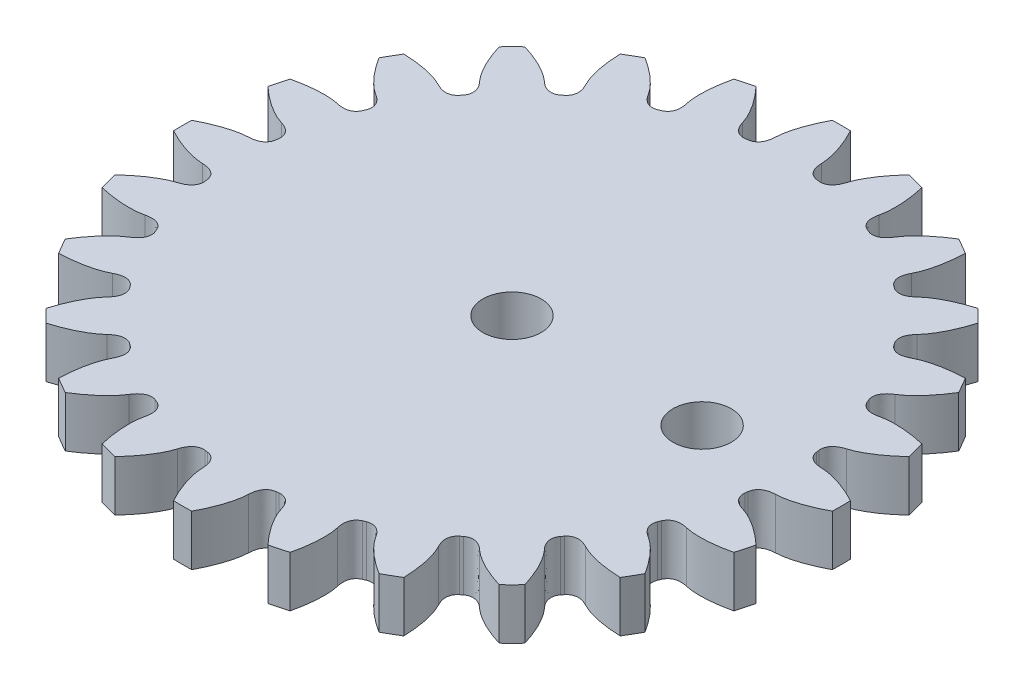
SolidWorks part; units mm, degrees
ref_plane "Спереди" through (0, 0, 0) normal (0, 0, 1) x (1, 0, 0)
ref_plane "Сверху" through (0, 0, 0) normal (0, 1, 0) x (1, 0, 0)
ref_plane "Справа" through (0, 0, 0) normal (1, 0, 0) x (0, 0, -1)
sketch "Эскиз1" plane through (0, 0, 0) normal (0, 1, 0) x (1, 0, 0)
  line L0 (0, 0) -> (7.5, 0) construction
  circle A0 centre (0, 0) radius 1.15
  circle A2 centre (7.5, 0) radius 1.15
  line B0 (-14.3, 0) -> (14.3, 0) construction
  line B1 (0, -14.3) -> (0, 14.3) construction
  arc B2 (0.3577, 12.9951) -> (-0.3577, 12.9951) centre (0, 0) ccw
  arc B3 (-1.346, 10.6654) -> (-1.4603, 10.6504) centre (0, 0) ccw
  arc B4 (-3.0178, 12.6449) -> (-3.7089, 12.4597) centre (0, 0) ccw
  arc B5 (-4.0605, 9.9536) -> (-4.1671, 9.9095) centre (0, 0) ccw
  arc B6 (-6.1877, 11.4329) -> (-6.8073, 11.0752) centre (0, 0) ccw
  arc B7 (-6.4984, 8.5635) -> (-6.5898, 8.4933) centre (0, 0) ccw
  arc B8 (-8.936, 9.4419) -> (-9.4419, 8.936) centre (0, 0) ccw
  arc B9 (-8.4933, 6.5898) -> (-8.5635, 6.4984) centre (0, 0) ccw
  arc B10 (-11.0752, 6.8073) -> (-11.4329, 6.1877) centre (0, 0) ccw
  arc B11 (-9.9095, 4.1671) -> (-9.9536, 4.0605) centre (0, 0) ccw
  arc B12 (-12.4597, 3.7089) -> (-12.6449, 3.0178) centre (0, 0) ccw
  arc B13 (-10.6504, 1.4603) -> (-10.6654, 1.346) centre (0, 0) ccw
  arc B14 (-12.9951, 0.3577) -> (-12.9951, -0.3577) centre (0, 0) ccw
  arc B15 (-10.6654, -1.346) -> (-10.6504, -1.4603) centre (0, 0) ccw
  arc B16 (-12.6449, -3.0178) -> (-12.4597, -3.7089) centre (0, 0) ccw
  arc B17 (-9.9536, -4.0605) -> (-9.9095, -4.1671) centre (0, 0) ccw
  arc B18 (-11.4329, -6.1877) -> (-11.0752, -6.8073) centre (0, 0) ccw
  arc B19 (-8.5635, -6.4984) -> (-8.4933, -6.5898) centre (0, 0) ccw
  arc B20 (-9.4419, -8.936) -> (-8.936, -9.4419) centre (0, 0) ccw
  arc B21 (-6.5898, -8.4933) -> (-6.4984, -8.5635) centre (0, 0) ccw
  arc B22 (-6.8073, -11.0752) -> (-6.1877, -11.4329) centre (0, 0) ccw
  arc B23 (-4.1671, -9.9095) -> (-4.0605, -9.9536) centre (0, 0) ccw
  arc B24 (-3.7089, -12.4597) -> (-3.0178, -12.6449) centre (0, 0) ccw
  arc B25 (-1.4603, -10.6504) -> (-1.346, -10.6654) centre (0, 0) ccw
  arc B26 (-0.3577, -12.9951) -> (0.3577, -12.9951) centre (0, 0) ccw
  arc B27 (1.346, -10.6654) -> (1.4603, -10.6504) centre (0, 0) ccw
  arc B28 (3.0178, -12.6449) -> (3.7089, -12.4597) centre (0, 0) ccw
  arc B29 (4.0605, -9.9536) -> (4.1671, -9.9095) centre (0, 0) ccw
  arc B30 (6.1877, -11.4329) -> (6.8073, -11.0752) centre (0, 0) ccw
  arc B31 (6.4984, -8.5635) -> (6.5898, -8.4933) centre (0, 0) ccw
  arc B32 (8.936, -9.4419) -> (9.4419, -8.936) centre (0, 0) ccw
  arc B33 (8.4933, -6.5898) -> (8.5635, -6.4984) centre (0, 0) ccw
  arc B34 (11.0752, -6.8073) -> (11.4329, -6.1877) centre (0, 0) ccw
  arc B35 (9.9095, -4.1671) -> (9.9536, -4.0605) centre (0, 0) ccw
  arc B36 (12.4597, -3.7089) -> (12.6449, -3.0178) centre (0, 0) ccw
  arc B37 (10.6504, -1.4603) -> (10.6654, -1.346) centre (0, 0) ccw
  arc B38 (12.9951, -0.3577) -> (12.9951, 0.3577) centre (0, 0) ccw
  arc B39 (10.6654, 1.346) -> (10.6504, 1.4603) centre (0, 0) ccw
  arc B40 (12.6449, 3.0178) -> (12.4597, 3.7089) centre (0, 0) ccw
  arc B41 (9.9536, 4.0605) -> (9.9095, 4.1671) centre (0, 0) ccw
  arc B42 (11.4329, 6.1877) -> (11.0752, 6.8073) centre (0, 0) ccw
  arc B43 (8.5635, 6.4984) -> (8.4933, 6.5898) centre (0, 0) ccw
  arc B44 (9.4419, 8.936) -> (8.936, 9.4419) centre (0, 0) ccw
  arc B45 (6.5898, 8.4933) -> (6.4984, 8.5635) centre (0, 0) ccw
  arc B46 (6.8073, 11.0752) -> (6.1877, 11.4329) centre (0, 0) ccw
  arc B47 (4.1671, 9.9095) -> (4.0605, 9.9536) centre (0, 0) ccw
  arc B48 (3.7089, 12.4597) -> (3.0178, 12.6449) centre (0, 0) ccw
  arc B49 (1.4603, 10.6504) -> (1.346, 10.6654) centre (0, 0) ccw
  circle B50 centre (0, 0) radius 12 construction
  spline B51 degree 3 poles (0.9058, 11.3017) (0.9058, 11.2304) (0.9138, 11.1608) (0.9299, 11.0929) (0.9396, 11.0522) (0.9513, 11.0113) (0.9676, 10.9727) (0.9799, 10.9437) (0.994, 10.915) (1.0107, 10.8883) (1.0248, 10.8656) (1.0406, 10.8436) (1.058, 10.8234) (1.0738, 10.805) (1.091, 10.7875) (1.1093, 10.7717) (1.1266, 10.7569) (1.1451, 10.7431) (1.1643, 10.7309) (1.1829, 10.7192) (1.2025, 10.7087) (1.2225, 10.6998) (1.2421, 10.6911) (1.2626, 10.6838) (1.2833, 10.678) (1.3038, 10.6723) (1.3247, 10.6681) (1.346, 10.6654) knots 0 0 0 0 1 1 1 2 2 2 3 3 3 4 4 4 5 5 5 6 6 6 7 7 7 8 8 8 9 9 9 9
  spline B52 degree 3 poles (-0.9058, 11.3017) (-0.9058, 11.2304) (-0.9138, 11.1608) (-0.9299, 11.0929) (-0.9396, 11.0522) (-0.9513, 11.0113) (-0.9676, 10.9727) (-0.9799, 10.9437) (-0.994, 10.915) (-1.0107, 10.8883) (-1.0248, 10.8656) (-1.0406, 10.8436) (-1.058, 10.8234) (-1.0738, 10.805) (-1.091, 10.7875) (-1.1093, 10.7717) (-1.1266, 10.7569) (-1.1451, 10.7431) (-1.1643, 10.7309) (-1.1829, 10.7192) (-1.2025, 10.7087) (-1.2225, 10.6998) (-1.2421, 10.6911) (-1.2626, 10.6838) (-1.2833, 10.678) (-1.3038, 10.6723) (-1.3247, 10.6681) (-1.346, 10.6654) knots 0 0 0 0 1 1 1 2 2 2 3 3 3 4 4 4 5 5 5 6 6 6 7 7 7 8 8 8 9 9 9 9
  spline B53 degree 3 poles (0.9058, 11.3017) (0.9032, 11.3642) (0.898, 11.4263) (0.8903, 11.4882) (0.8824, 11.551) (0.8712, 11.6136) (0.8589, 11.6757) (0.8463, 11.7389) (0.8314, 11.8016) (0.8153, 11.864) (0.7989, 11.9273) (0.7806, 11.9902) (0.7612, 12.0526) (0.7414, 12.116) (0.72, 12.179) (0.6975, 12.2415) (0.6746, 12.3049) (0.6503, 12.3678) (0.6249, 12.4303) (0.5991, 12.4937) (0.572, 12.5566) (0.5439, 12.6189) (0.5153, 12.6822) (0.4855, 12.745) (0.4547, 12.8073) (0.4235, 12.8704) (0.3912, 12.933) (0.3577, 12.9951) knots 0 0 0 0 1 1 1 2 2 2 3 3 3 4 4 4 5 5 5 6 6 6 7 7 7 8 8 8 9 9 9 9
  spline B54 degree 3 poles (-0.9058, 11.3017) (-0.9032, 11.3642) (-0.898, 11.4263) (-0.8903, 11.4882) (-0.8824, 11.551) (-0.8712, 11.6136) (-0.8589, 11.6757) (-0.8463, 11.7389) (-0.8314, 11.8016) (-0.8153, 11.864) (-0.7989, 11.9273) (-0.7806, 11.9902) (-0.7612, 12.0526) (-0.7414, 12.116) (-0.72, 12.179) (-0.6975, 12.2415) (-0.6746, 12.3049) (-0.6503, 12.3678) (-0.6249, 12.4303) (-0.5991, 12.4937) (-0.572, 12.5566) (-0.5439, 12.6189) (-0.5153, 12.6822) (-0.4855, 12.745) (-0.4547, 12.8073) (-0.4235, 12.8704) (-0.3912, 12.933) (-0.3577, 12.9951) knots 0 0 0 0 1 1 1 2 2 2 3 3 3 4 4 4 5 5 5 6 6 6 7 7 7 8 8 8 9 9 9 9
  spline B55 degree 3 poles (-2.0502, 11.151) (-2.0317, 11.0822) (-2.0059, 11.017) (-1.9728, 10.9556) (-1.9529, 10.9188) (-1.931, 10.8823) (-1.9053, 10.8493) (-1.886, 10.8244) (-1.8649, 10.8004) (-1.8419, 10.7789) (-1.8224, 10.7606) (-1.8014, 10.7435) (-1.7793, 10.7284) (-1.7594, 10.7148) (-1.7382, 10.7023) (-1.7164, 10.6918) (-1.6959, 10.6819) (-1.6745, 10.6734) (-1.6527, 10.6666) (-1.6318, 10.6601) (-1.6101, 10.655) (-1.5885, 10.6516) (-1.5672, 10.6483) (-1.5456, 10.6465) (-1.5241, 10.6463) (-1.5028, 10.6461) (-1.4816, 10.6475) (-1.4603, 10.6504) knots 0 0 0 0 1 1 1 2 2 2 3 3 3 4 4 4 5 5 5 6 6 6 7 7 7 8 8 8 9 9 9 9
  spline B56 degree 3 poles (-3.8, 10.6822) (-3.7815, 10.6133) (-3.7713, 10.544) (-3.7693, 10.4743) (-3.7681, 10.4325) (-3.7688, 10.3898) (-3.7746, 10.3484) (-3.7789, 10.3172) (-3.7852, 10.2858) (-3.7943, 10.2557) (-3.8021, 10.2302) (-3.8117, 10.2048) (-3.8232, 10.1807) (-3.8337, 10.1589) (-3.8458, 10.1376) (-3.8595, 10.1176) (-3.8723, 10.0988) (-3.8866, 10.0806) (-3.902, 10.0639) (-3.9169, 10.0478) (-3.9331, 10.0326) (-3.9502, 10.0188) (-3.9669, 10.0053) (-3.9848, 9.9929) (-4.0032, 9.982) (-4.0216, 9.9712) (-4.0406, 9.9618) (-4.0605, 9.9536) knots 0 0 0 0 1 1 1 2 2 2 3 3 3 4 4 4 5 5 5 6 6 6 7 7 7 8 8 8 9 9 9 9
  spline B57 degree 3 poles (-2.0502, 11.151) (-2.0689, 11.2107) (-2.09, 11.2694) (-2.1134, 11.3271) (-2.1373, 11.3858) (-2.1643, 11.4434) (-2.1923, 11.5002) (-2.2208, 11.5579) (-2.2514, 11.6147) (-2.2831, 11.6707) (-2.3153, 11.7276) (-2.3493, 11.7837) (-2.3842, 11.8389) (-2.4197, 11.8951) (-2.4567, 11.9503) (-2.4946, 12.0049) (-2.5331, 12.0602) (-2.5729, 12.1147) (-2.6136, 12.1685) (-2.6549, 12.223) (-2.6974, 12.2768) (-2.7407, 12.3297) (-2.7847, 12.3835) (-2.8297, 12.4364) (-2.8755, 12.4885) (-2.9221, 12.5415) (-2.9695, 12.5936) (-3.0178, 12.6449) knots 0 0 0 0 1 1 1 2 2 2 3 3 3 4 4 4 5 5 5 6 6 6 7 7 7 8 8 8 9 9 9 9
  spline B58 degree 3 poles (-3.8, 10.6822) (-3.8136, 10.7432) (-3.8247, 10.8046) (-3.8333, 10.8663) (-3.842, 10.929) (-3.8474, 10.9924) (-3.8515, 11.0556) (-3.8557, 11.1198) (-3.8576, 11.1843) (-3.8581, 11.2487) (-3.8587, 11.3141) (-3.8573, 11.3796) (-3.8547, 11.4449) (-3.852, 11.5113) (-3.8476, 11.5776) (-3.8421, 11.6438) (-3.8364, 11.711) (-3.8292, 11.7781) (-3.8208, 11.845) (-3.8123, 11.9129) (-3.8024, 11.9807) (-3.7914, 12.0482) (-3.7802, 12.1167) (-3.7676, 12.1851) (-3.754, 12.2532) (-3.7402, 12.3223) (-3.7251, 12.3911) (-3.7089, 12.4597) knots 0 0 0 0 1 1 1 2 2 2 3 3 3 4 4 4 5 5 5 6 6 6 7 7 7 8 8 8 9 9 9 9
  spline B59 degree 3 poles (-4.8664, 10.2404) (-4.8308, 10.1787) (-4.789, 10.1225) (-4.7411, 10.0717) (-4.7124, 10.0413) (-4.6817, 10.0117) (-4.6484, 9.9865) (-4.6233, 9.9675) (-4.5967, 9.9497) (-4.5689, 9.9349) (-4.5453, 9.9223) (-4.5206, 9.9111) (-4.4954, 9.9023) (-4.4726, 9.8943) (-4.4489, 9.8878) (-4.4252, 9.8833) (-4.4028, 9.879) (-4.3799, 9.8763) (-4.3571, 9.8754) (-4.3352, 9.8745) (-4.313, 9.8752) (-4.2912, 9.8776) (-4.2698, 9.8798) (-4.2484, 9.8837) (-4.2276, 9.8891) (-4.2071, 9.8944) (-4.1869, 9.9012) (-4.1671, 9.9095) knots 0 0 0 0 1 1 1 2 2 2 3 3 3 4 4 4 5 5 5 6 6 6 7 7 7 8 8 8 9 9 9 9
  spline B60 degree 3 poles (-6.4353, 9.3347) (-6.3996, 9.2729) (-6.3718, 9.2086) (-6.3518, 9.1418) (-6.3398, 9.1017) (-6.3295, 9.0604) (-6.3243, 9.0188) (-6.3204, 8.9876) (-6.3184, 8.9557) (-6.3194, 8.9242) (-6.3203, 8.8975) (-6.323, 8.8706) (-6.3279, 8.8443) (-6.3324, 8.8205) (-6.3386, 8.7968) (-6.3466, 8.7739) (-6.3541, 8.7524) (-6.3632, 8.7312) (-6.3738, 8.7111) (-6.384, 8.6917) (-6.3957, 8.6728) (-6.4086, 8.655) (-6.4213, 8.6377) (-6.4353, 8.6211) (-6.4504, 8.6058) (-6.4653, 8.5906) (-6.4813, 8.5765) (-6.4984, 8.5635) knots 0 0 0 0 1 1 1 2 2 2 3 3 3 4 4 4 5 5 5 6 6 6 7 7 7 8 8 8 9 9 9 9
  spline B61 degree 3 poles (-4.8664, 10.2404) (-4.8999, 10.2932) (-4.9355, 10.3445) (-4.9731, 10.3942) (-5.0113, 10.4447) (-5.0523, 10.4933) (-5.0941, 10.5409) (-5.1365, 10.5893) (-5.1808, 10.6362) (-5.2259, 10.6822) (-5.2718, 10.7288) (-5.319, 10.7741) (-5.3671, 10.8185) (-5.4159, 10.8635) (-5.4659, 10.9073) (-5.5167, 10.9502) (-5.5682, 10.9937) (-5.6207, 11.036) (-5.674, 11.0774) (-5.728, 11.1194) (-5.7829, 11.1603) (-5.8385, 11.2003) (-5.8949, 11.2408) (-5.9521, 11.2803) (-6.0098, 11.3188) (-6.0685, 11.3578) (-6.1278, 11.3959) (-6.1877, 11.4329) knots 0 0 0 0 1 1 1 2 2 2 3 3 3 4 4 4 5 5 5 6 6 6 7 7 7 8 8 8 9 9 9 9
  spline B62 degree 3 poles (-6.4353, 9.3347) (-6.4642, 9.3901) (-6.4908, 9.4465) (-6.5151, 9.5039) (-6.5397, 9.5623) (-6.5613, 9.622) (-6.5817, 9.6821) (-6.6024, 9.743) (-6.6209, 9.8048) (-6.638, 9.8669) (-6.6555, 9.9299) (-6.6711, 9.9935) (-6.6855, 10.0573) (-6.7001, 10.1221) (-6.713, 10.1873) (-6.7248, 10.2527) (-6.7367, 10.319) (-6.7471, 10.3857) (-6.7563, 10.4525) (-6.7657, 10.5203) (-6.7737, 10.5883) (-6.7805, 10.6564) (-6.7874, 10.7255) (-6.793, 10.7948) (-6.7974, 10.8641) (-6.8019, 10.9344) (-6.8053, 11.0047) (-6.8073, 11.0752) knots 0 0 0 0 1 1 1 2 2 2 3 3 3 4 4 4 5 5 5 6 6 6 7 7 7 8 8 8 9 9 9 9
  spline B63 degree 3 poles (-7.351, 8.632) (-7.3006, 8.5816) (-7.2457, 8.5381) (-7.1863, 8.5015) (-7.1507, 8.4795) (-7.1134, 8.4588) (-7.0747, 8.4431) (-7.0455, 8.4312) (-7.0152, 8.421) (-6.9845, 8.4138) (-6.9585, 8.4078) (-6.9318, 8.4034) (-6.9052, 8.4014) (-6.881, 8.3996) (-6.8565, 8.3994) (-6.8324, 8.4012) (-6.8097, 8.4029) (-6.7868, 8.4062) (-6.7646, 8.4112) (-6.7432, 8.416) (-6.7219, 8.4224) (-6.7015, 8.4304) (-6.6814, 8.4381) (-6.6618, 8.4474) (-6.6431, 8.4579) (-6.6246, 8.4684) (-6.6068, 8.4802) (-6.5898, 8.4933) knots 0 0 0 0 1 1 1 2 2 2 3 3 3 4 4 4 5 5 5 6 6 6 7 7 7 8 8 8 9 9 9 9
  spline B64 degree 3 poles (-8.632, 7.351) (-8.5816, 7.3006) (-8.5381, 7.2457) (-8.5015, 7.1863) (-8.4795, 7.1507) (-8.4588, 7.1134) (-8.4431, 7.0747) (-8.4312, 7.0455) (-8.421, 7.0152) (-8.4138, 6.9845) (-8.4078, 6.9585) (-8.4034, 6.9318) (-8.4014, 6.9052) (-8.3996, 6.881) (-8.3994, 6.8565) (-8.4012, 6.8324) (-8.4029, 6.8097) (-8.4062, 6.7868) (-8.4112, 6.7646) (-8.416, 6.7432) (-8.4224, 6.7219) (-8.4304, 6.7015) (-8.4381, 6.6814) (-8.4474, 6.6618) (-8.4579, 6.6431) (-8.4684, 6.6246) (-8.4802, 6.6068) (-8.4933, 6.5898) knots 0 0 0 0 1 1 1 2 2 2 3 3 3 4 4 4 5 5 5 6 6 6 7 7 7 8 8 8 9 9 9 9
  spline B65 degree 3 poles (-7.351, 8.632) (-7.3971, 8.6743) (-7.4447, 8.7146) (-7.4938, 8.7529) (-7.5438, 8.7918) (-7.596, 8.8281) (-7.6487, 8.8633) (-7.7022, 8.8991) (-7.7571, 8.9329) (-7.8126, 8.9656) (-7.869, 8.9988) (-7.9263, 9.0303) (-7.9843, 9.0607) (-8.0431, 9.0916) (-8.1027, 9.121) (-8.1628, 9.1492) (-8.2238, 9.1779) (-8.2855, 9.2052) (-8.3477, 9.2314) (-8.4107, 9.258) (-8.4744, 9.2833) (-8.5384, 9.3075) (-8.6033, 9.3321) (-8.6688, 9.3554) (-8.7346, 9.3776) (-8.8013, 9.4002) (-8.8684, 9.4216) (-8.936, 9.4419) knots 0 0 0 0 1 1 1 2 2 2 3 3 3 4 4 4 5 5 5 6 6 6 7 7 7 8 8 8 9 9 9 9
  spline B66 degree 3 poles (-8.632, 7.351) (-8.6743, 7.3971) (-8.7146, 7.4447) (-8.7529, 7.4938) (-8.7918, 7.5438) (-8.8281, 7.596) (-8.8633, 7.6487) (-8.8991, 7.7022) (-8.9329, 7.7571) (-8.9656, 7.8126) (-8.9988, 7.869) (-9.0303, 7.9263) (-9.0607, 7.9843) (-9.0916, 8.0431) (-9.121, 8.1027) (-9.1492, 8.1628) (-9.1779, 8.2238) (-9.2052, 8.2855) (-9.2314, 8.3477) (-9.258, 8.4107) (-9.2833, 8.4744) (-9.3075, 8.5384) (-9.3321, 8.6033) (-9.3554, 8.6688) (-9.3776, 8.7346) (-9.4002, 8.8013) (-9.4216, 8.8684) (-9.4419, 8.936) knots 0 0 0 0 1 1 1 2 2 2 3 3 3 4 4 4 5 5 5 6 6 6 7 7 7 8 8 8 9 9 9 9
  spline B67 degree 3 poles (-9.3347, 6.4353) (-9.2729, 6.3996) (-9.2086, 6.3718) (-9.1418, 6.3518) (-9.1017, 6.3398) (-9.0604, 6.3295) (-9.0188, 6.3243) (-8.9876, 6.3204) (-8.9557, 6.3184) (-8.9242, 6.3194) (-8.8975, 6.3203) (-8.8706, 6.323) (-8.8443, 6.3279) (-8.8205, 6.3324) (-8.7968, 6.3386) (-8.7739, 6.3466) (-8.7524, 6.3541) (-8.7312, 6.3632) (-8.7111, 6.3738) (-8.6917, 6.384) (-8.6728, 6.3957) (-8.655, 6.4086) (-8.6377, 6.4213) (-8.6211, 6.4353) (-8.6058, 6.4504) (-8.5906, 6.4653) (-8.5765, 6.4813) (-8.5635, 6.4984) knots 0 0 0 0 1 1 1 2 2 2 3 3 3 4 4 4 5 5 5 6 6 6 7 7 7 8 8 8 9 9 9 9
  spline B68 degree 3 poles (-10.2404, 4.8664) (-10.1787, 4.8308) (-10.1225, 4.789) (-10.0717, 4.7411) (-10.0413, 4.7124) (-10.0117, 4.6817) (-9.9865, 4.6484) (-9.9675, 4.6233) (-9.9497, 4.5967) (-9.9349, 4.5689) (-9.9223, 4.5453) (-9.9111, 4.5206) (-9.9023, 4.4954) (-9.8943, 4.4726) (-9.8878, 4.4489) (-9.8833, 4.4252) (-9.879, 4.4028) (-9.8763, 4.3799) (-9.8754, 4.3571) (-9.8745, 4.3352) (-9.8752, 4.313) (-9.8776, 4.2912) (-9.8798, 4.2698) (-9.8837, 4.2484) (-9.8891, 4.2276) (-9.8944, 4.2071) (-9.9012, 4.1869) (-9.9095, 4.1671) knots 0 0 0 0 1 1 1 2 2 2 3 3 3 4 4 4 5 5 5 6 6 6 7 7 7 8 8 8 9 9 9 9
  spline B69 degree 3 poles (-9.3347, 6.4353) (-9.3901, 6.4642) (-9.4465, 6.4908) (-9.5039, 6.5151) (-9.5623, 6.5397) (-9.622, 6.5613) (-9.6821, 6.5817) (-9.743, 6.6024) (-9.8048, 6.6209) (-9.8669, 6.638) (-9.9299, 6.6555) (-9.9935, 6.6711) (-10.0573, 6.6855) (-10.1221, 6.7001) (-10.1873, 6.713) (-10.2527, 6.7248) (-10.319, 6.7367) (-10.3857, 6.7471) (-10.4525, 6.7563) (-10.5203, 6.7657) (-10.5883, 6.7737) (-10.6564, 6.7805) (-10.7255, 6.7874) (-10.7948, 6.793) (-10.8641, 6.7974) (-10.9344, 6.8019) (-11.0047, 6.8053) (-11.0752, 6.8073) knots 0 0 0 0 1 1 1 2 2 2 3 3 3 4 4 4 5 5 5 6 6 6 7 7 7 8 8 8 9 9 9 9
  spline B70 degree 3 poles (-10.2404, 4.8664) (-10.2932, 4.8999) (-10.3445, 4.9355) (-10.3942, 4.9731) (-10.4447, 5.0113) (-10.4933, 5.0523) (-10.5409, 5.0941) (-10.5893, 5.1365) (-10.6362, 5.1808) (-10.6822, 5.2259) (-10.7288, 5.2718) (-10.7741, 5.319) (-10.8185, 5.3671) (-10.8635, 5.4159) (-10.9073, 5.4659) (-10.9502, 5.5167) (-10.9937, 5.5682) (-11.036, 5.6207) (-11.0774, 5.674) (-11.1194, 5.728) (-11.1603, 5.7829) (-11.2003, 5.8385) (-11.2408, 5.8949) (-11.2803, 5.9521) (-11.3188, 6.0098) (-11.3578, 6.0685) (-11.3959, 6.1278) (-11.4329, 6.1877) knots 0 0 0 0 1 1 1 2 2 2 3 3 3 4 4 4 5 5 5 6 6 6 7 7 7 8 8 8 9 9 9 9
  spline B71 degree 3 poles (-10.6822, 3.8) (-10.6133, 3.7815) (-10.544, 3.7713) (-10.4743, 3.7693) (-10.4325, 3.7681) (-10.3898, 3.7688) (-10.3484, 3.7746) (-10.3172, 3.7789) (-10.2858, 3.7852) (-10.2557, 3.7943) (-10.2302, 3.8021) (-10.2048, 3.8117) (-10.1807, 3.8232) (-10.1589, 3.8337) (-10.1376, 3.8458) (-10.1176, 3.8595) (-10.0988, 3.8723) (-10.0806, 3.8866) (-10.0639, 3.902) (-10.0478, 3.9169) (-10.0326, 3.9331) (-10.0188, 3.9502) (-10.0053, 3.9669) (-9.9929, 3.9848) (-9.982, 4.0032) (-9.9712, 4.0216) (-9.9618, 4.0406) (-9.9536, 4.0605) knots 0 0 0 0 1 1 1 2 2 2 3 3 3 4 4 4 5 5 5 6 6 6 7 7 7 8 8 8 9 9 9 9
  spline B72 degree 3 poles (-11.151, 2.0502) (-11.0822, 2.0317) (-11.017, 2.0059) (-10.9556, 1.9728) (-10.9188, 1.9529) (-10.8823, 1.931) (-10.8493, 1.9053) (-10.8244, 1.886) (-10.8004, 1.8649) (-10.7789, 1.8419) (-10.7606, 1.8224) (-10.7435, 1.8014) (-10.7284, 1.7793) (-10.7148, 1.7594) (-10.7023, 1.7382) (-10.6918, 1.7164) (-10.6819, 1.6959) (-10.6734, 1.6745) (-10.6666, 1.6527) (-10.6601, 1.6318) (-10.655, 1.6101) (-10.6516, 1.5885) (-10.6483, 1.5672) (-10.6465, 1.5456) (-10.6463, 1.5241) (-10.6461, 1.5028) (-10.6475, 1.4816) (-10.6504, 1.4603) knots 0 0 0 0 1 1 1 2 2 2 3 3 3 4 4 4 5 5 5 6 6 6 7 7 7 8 8 8 9 9 9 9
  spline B73 degree 3 poles (-10.6822, 3.8) (-10.7432, 3.8136) (-10.8046, 3.8247) (-10.8663, 3.8333) (-10.929, 3.842) (-10.9924, 3.8474) (-11.0556, 3.8515) (-11.1198, 3.8557) (-11.1843, 3.8576) (-11.2487, 3.8581) (-11.3141, 3.8587) (-11.3796, 3.8573) (-11.4449, 3.8547) (-11.5113, 3.852) (-11.5776, 3.8476) (-11.6438, 3.8421) (-11.711, 3.8364) (-11.7781, 3.8292) (-11.845, 3.8208) (-11.9129, 3.8123) (-11.9807, 3.8024) (-12.0482, 3.7914) (-12.1167, 3.7802) (-12.1851, 3.7676) (-12.2532, 3.754) (-12.3223, 3.7402) (-12.3911, 3.7251) (-12.4597, 3.7089) knots 0 0 0 0 1 1 1 2 2 2 3 3 3 4 4 4 5 5 5 6 6 6 7 7 7 8 8 8 9 9 9 9
  spline B74 degree 3 poles (-11.151, 2.0502) (-11.2107, 2.0689) (-11.2694, 2.09) (-11.3271, 2.1134) (-11.3858, 2.1373) (-11.4434, 2.1643) (-11.5002, 2.1923) (-11.5579, 2.2208) (-11.6147, 2.2514) (-11.6707, 2.2831) (-11.7276, 2.3153) (-11.7837, 2.3493) (-11.8389, 2.3842) (-11.8951, 2.4197) (-11.9503, 2.4567) (-12.0049, 2.4946) (-12.0602, 2.5331) (-12.1147, 2.5729) (-12.1685, 2.6136) (-12.223, 2.6549) (-12.2768, 2.6974) (-12.3297, 2.7407) (-12.3835, 2.7847) (-12.4364, 2.8297) (-12.4885, 2.8755) (-12.5415, 2.9221) (-12.5936, 2.9695) (-12.6449, 3.0178) knots 0 0 0 0 1 1 1 2 2 2 3 3 3 4 4 4 5 5 5 6 6 6 7 7 7 8 8 8 9 9 9 9
  spline B75 degree 3 poles (-11.3017, 0.9058) (-11.2304, 0.9058) (-11.1608, 0.9138) (-11.0929, 0.9299) (-11.0522, 0.9396) (-11.0113, 0.9513) (-10.9727, 0.9676) (-10.9437, 0.9799) (-10.915, 0.994) (-10.8883, 1.0107) (-10.8656, 1.0248) (-10.8436, 1.0406) (-10.8234, 1.058) (-10.805, 1.0738) (-10.7875, 1.091) (-10.7717, 1.1093) (-10.7569, 1.1266) (-10.7431, 1.1451) (-10.7309, 1.1643) (-10.7192, 1.1829) (-10.7087, 1.2025) (-10.6998, 1.2225) (-10.6911, 1.2421) (-10.6838, 1.2626) (-10.678, 1.2833) (-10.6723, 1.3038) (-10.6681, 1.3247) (-10.6654, 1.346) knots 0 0 0 0 1 1 1 2 2 2 3 3 3 4 4 4 5 5 5 6 6 6 7 7 7 8 8 8 9 9 9 9
  spline B76 degree 3 poles (-11.3017, -0.9058) (-11.2304, -0.9058) (-11.1608, -0.9138) (-11.0929, -0.9299) (-11.0522, -0.9396) (-11.0113, -0.9513) (-10.9727, -0.9676) (-10.9437, -0.9799) (-10.915, -0.994) (-10.8883, -1.0107) (-10.8656, -1.0248) (-10.8436, -1.0406) (-10.8234, -1.058) (-10.805, -1.0738) (-10.7875, -1.091) (-10.7717, -1.1093) (-10.7569, -1.1266) (-10.7431, -1.1451) (-10.7309, -1.1643) (-10.7192, -1.1829) (-10.7087, -1.2025) (-10.6998, -1.2225) (-10.6911, -1.2421) (-10.6838, -1.2626) (-10.678, -1.2833) (-10.6723, -1.3038) (-10.6681, -1.3247) (-10.6654, -1.346) knots 0 0 0 0 1 1 1 2 2 2 3 3 3 4 4 4 5 5 5 6 6 6 7 7 7 8 8 8 9 9 9 9
  spline B77 degree 3 poles (-11.3017, 0.9058) (-11.3642, 0.9032) (-11.4263, 0.898) (-11.4882, 0.8903) (-11.551, 0.8824) (-11.6136, 0.8712) (-11.6757, 0.8589) (-11.7389, 0.8463) (-11.8016, 0.8314) (-11.864, 0.8153) (-11.9273, 0.7989) (-11.9902, 0.7806) (-12.0526, 0.7612) (-12.116, 0.7414) (-12.179, 0.72) (-12.2415, 0.6975) (-12.3049, 0.6746) (-12.3678, 0.6503) (-12.4303, 0.6249) (-12.4937, 0.5991) (-12.5566, 0.572) (-12.6189, 0.5439) (-12.6822, 0.5153) (-12.745, 0.4855) (-12.8073, 0.4547) (-12.8704, 0.4235) (-12.933, 0.3912) (-12.9951, 0.3577) knots 0 0 0 0 1 1 1 2 2 2 3 3 3 4 4 4 5 5 5 6 6 6 7 7 7 8 8 8 9 9 9 9
  spline B78 degree 3 poles (-11.3017, -0.9058) (-11.3642, -0.9032) (-11.4263, -0.898) (-11.4882, -0.8903) (-11.551, -0.8824) (-11.6136, -0.8712) (-11.6757, -0.8589) (-11.7389, -0.8463) (-11.8016, -0.8314) (-11.864, -0.8153) (-11.9273, -0.7989) (-11.9902, -0.7806) (-12.0526, -0.7612) (-12.116, -0.7414) (-12.179, -0.72) (-12.2415, -0.6975) (-12.3049, -0.6746) (-12.3678, -0.6503) (-12.4303, -0.6249) (-12.4937, -0.5991) (-12.5566, -0.572) (-12.6189, -0.5439) (-12.6822, -0.5153) (-12.745, -0.4855) (-12.8073, -0.4547) (-12.8704, -0.4235) (-12.933, -0.3912) (-12.9951, -0.3577) knots 0 0 0 0 1 1 1 2 2 2 3 3 3 4 4 4 5 5 5 6 6 6 7 7 7 8 8 8 9 9 9 9
  spline B79 degree 3 poles (-11.151, -2.0502) (-11.0822, -2.0317) (-11.017, -2.0059) (-10.9556, -1.9728) (-10.9188, -1.9529) (-10.8823, -1.931) (-10.8493, -1.9053) (-10.8244, -1.886) (-10.8004, -1.8649) (-10.7789, -1.8419) (-10.7606, -1.8224) (-10.7435, -1.8014) (-10.7284, -1.7793) (-10.7148, -1.7594) (-10.7023, -1.7382) (-10.6918, -1.7164) (-10.6819, -1.6959) (-10.6734, -1.6745) (-10.6666, -1.6527) (-10.6601, -1.6318) (-10.655, -1.6101) (-10.6516, -1.5885) (-10.6483, -1.5672) (-10.6465, -1.5456) (-10.6463, -1.5241) (-10.6461, -1.5028) (-10.6475, -1.4816) (-10.6504, -1.4603) knots 0 0 0 0 1 1 1 2 2 2 3 3 3 4 4 4 5 5 5 6 6 6 7 7 7 8 8 8 9 9 9 9
  spline B80 degree 3 poles (-10.6822, -3.8) (-10.6133, -3.7815) (-10.544, -3.7713) (-10.4743, -3.7693) (-10.4325, -3.7681) (-10.3898, -3.7688) (-10.3484, -3.7746) (-10.3172, -3.7789) (-10.2858, -3.7852) (-10.2557, -3.7943) (-10.2302, -3.8021) (-10.2048, -3.8117) (-10.1807, -3.8232) (-10.1589, -3.8337) (-10.1376, -3.8458) (-10.1176, -3.8595) (-10.0988, -3.8723) (-10.0806, -3.8866) (-10.0639, -3.902) (-10.0478, -3.9169) (-10.0326, -3.9331) (-10.0188, -3.9502) (-10.0053, -3.9669) (-9.9929, -3.9848) (-9.982, -4.0032) (-9.9712, -4.0216) (-9.9618, -4.0406) (-9.9536, -4.0605) knots 0 0 0 0 1 1 1 2 2 2 3 3 3 4 4 4 5 5 5 6 6 6 7 7 7 8 8 8 9 9 9 9
  spline B81 degree 3 poles (-11.151, -2.0502) (-11.2107, -2.0689) (-11.2694, -2.09) (-11.3271, -2.1134) (-11.3858, -2.1373) (-11.4434, -2.1643) (-11.5002, -2.1923) (-11.5579, -2.2208) (-11.6147, -2.2514) (-11.6707, -2.2831) (-11.7276, -2.3153) (-11.7837, -2.3493) (-11.8389, -2.3842) (-11.8951, -2.4197) (-11.9503, -2.4567) (-12.0049, -2.4946) (-12.0602, -2.5331) (-12.1147, -2.5729) (-12.1685, -2.6136) (-12.223, -2.6549) (-12.2768, -2.6974) (-12.3297, -2.7407) (-12.3835, -2.7847) (-12.4364, -2.8297) (-12.4885, -2.8755) (-12.5415, -2.9221) (-12.5936, -2.9695) (-12.6449, -3.0178) knots 0 0 0 0 1 1 1 2 2 2 3 3 3 4 4 4 5 5 5 6 6 6 7 7 7 8 8 8 9 9 9 9
  spline B82 degree 3 poles (-10.6822, -3.8) (-10.7432, -3.8136) (-10.8046, -3.8247) (-10.8663, -3.8333) (-10.929, -3.842) (-10.9924, -3.8474) (-11.0556, -3.8515) (-11.1198, -3.8557) (-11.1843, -3.8576) (-11.2487, -3.8581) (-11.3141, -3.8587) (-11.3796, -3.8573) (-11.4449, -3.8547) (-11.5113, -3.852) (-11.5776, -3.8476) (-11.6438, -3.8421) (-11.711, -3.8364) (-11.7781, -3.8292) (-11.845, -3.8208) (-11.9129, -3.8123) (-11.9807, -3.8024) (-12.0482, -3.7914) (-12.1167, -3.7802) (-12.1851, -3.7676) (-12.2532, -3.754) (-12.3223, -3.7402) (-12.3911, -3.7251) (-12.4597, -3.7089) knots 0 0 0 0 1 1 1 2 2 2 3 3 3 4 4 4 5 5 5 6 6 6 7 7 7 8 8 8 9 9 9 9
  spline B83 degree 3 poles (-10.2404, -4.8664) (-10.1787, -4.8308) (-10.1225, -4.789) (-10.0717, -4.7411) (-10.0413, -4.7124) (-10.0117, -4.6817) (-9.9865, -4.6484) (-9.9675, -4.6233) (-9.9497, -4.5967) (-9.9349, -4.5689) (-9.9223, -4.5453) (-9.9111, -4.5206) (-9.9023, -4.4954) (-9.8943, -4.4726) (-9.8878, -4.4489) (-9.8833, -4.4252) (-9.879, -4.4028) (-9.8763, -4.3799) (-9.8754, -4.3571) (-9.8745, -4.3352) (-9.8752, -4.313) (-9.8776, -4.2912) (-9.8798, -4.2698) (-9.8837, -4.2484) (-9.8891, -4.2276) (-9.8944, -4.2071) (-9.9012, -4.1869) (-9.9095, -4.1671) knots 0 0 0 0 1 1 1 2 2 2 3 3 3 4 4 4 5 5 5 6 6 6 7 7 7 8 8 8 9 9 9 9
  spline B84 degree 3 poles (-9.3347, -6.4353) (-9.2729, -6.3996) (-9.2086, -6.3718) (-9.1418, -6.3518) (-9.1017, -6.3398) (-9.0604, -6.3295) (-9.0188, -6.3243) (-8.9876, -6.3204) (-8.9557, -6.3184) (-8.9242, -6.3194) (-8.8975, -6.3203) (-8.8706, -6.323) (-8.8443, -6.3279) (-8.8205, -6.3324) (-8.7968, -6.3386) (-8.7739, -6.3466) (-8.7524, -6.3541) (-8.7312, -6.3632) (-8.7111, -6.3738) (-8.6917, -6.384) (-8.6728, -6.3957) (-8.655, -6.4086) (-8.6377, -6.4213) (-8.6211, -6.4353) (-8.6058, -6.4504) (-8.5906, -6.4653) (-8.5765, -6.4813) (-8.5635, -6.4984) knots 0 0 0 0 1 1 1 2 2 2 3 3 3 4 4 4 5 5 5 6 6 6 7 7 7 8 8 8 9 9 9 9
  spline B85 degree 3 poles (-10.2404, -4.8664) (-10.2932, -4.8999) (-10.3445, -4.9355) (-10.3942, -4.9731) (-10.4447, -5.0113) (-10.4933, -5.0523) (-10.5409, -5.0941) (-10.5893, -5.1365) (-10.6362, -5.1808) (-10.6822, -5.2259) (-10.7288, -5.2718) (-10.7741, -5.319) (-10.8185, -5.3671) (-10.8635, -5.4159) (-10.9073, -5.4659) (-10.9502, -5.5167) (-10.9937, -5.5682) (-11.036, -5.6207) (-11.0774, -5.674) (-11.1194, -5.728) (-11.1603, -5.7829) (-11.2003, -5.8385) (-11.2408, -5.8949) (-11.2803, -5.9521) (-11.3188, -6.0098) (-11.3578, -6.0685) (-11.3959, -6.1278) (-11.4329, -6.1877) knots 0 0 0 0 1 1 1 2 2 2 3 3 3 4 4 4 5 5 5 6 6 6 7 7 7 8 8 8 9 9 9 9
  spline B86 degree 3 poles (-9.3347, -6.4353) (-9.3901, -6.4642) (-9.4465, -6.4908) (-9.5039, -6.5151) (-9.5623, -6.5397) (-9.622, -6.5613) (-9.6821, -6.5817) (-9.743, -6.6024) (-9.8048, -6.6209) (-9.8669, -6.638) (-9.9299, -6.6555) (-9.9935, -6.6711) (-10.0573, -6.6855) (-10.1221, -6.7001) (-10.1873, -6.713) (-10.2527, -6.7248) (-10.319, -6.7367) (-10.3857, -6.7471) (-10.4525, -6.7563) (-10.5203, -6.7657) (-10.5883, -6.7737) (-10.6564, -6.7805) (-10.7255, -6.7874) (-10.7948, -6.793) (-10.8641, -6.7974) (-10.9344, -6.8019) (-11.0047, -6.8053) (-11.0752, -6.8073) knots 0 0 0 0 1 1 1 2 2 2 3 3 3 4 4 4 5 5 5 6 6 6 7 7 7 8 8 8 9 9 9 9
  spline B87 degree 3 poles (-8.632, -7.351) (-8.5816, -7.3006) (-8.5381, -7.2457) (-8.5015, -7.1863) (-8.4795, -7.1507) (-8.4588, -7.1134) (-8.4431, -7.0747) (-8.4312, -7.0455) (-8.421, -7.0152) (-8.4138, -6.9845) (-8.4078, -6.9585) (-8.4034, -6.9318) (-8.4014, -6.9052) (-8.3996, -6.881) (-8.3994, -6.8565) (-8.4012, -6.8324) (-8.4029, -6.8097) (-8.4062, -6.7868) (-8.4112, -6.7646) (-8.416, -6.7432) (-8.4224, -6.7219) (-8.4304, -6.7015) (-8.4381, -6.6814) (-8.4474, -6.6618) (-8.4579, -6.6431) (-8.4684, -6.6246) (-8.4802, -6.6068) (-8.4933, -6.5898) knots 0 0 0 0 1 1 1 2 2 2 3 3 3 4 4 4 5 5 5 6 6 6 7 7 7 8 8 8 9 9 9 9
  spline B88 degree 3 poles (-7.351, -8.632) (-7.3006, -8.5816) (-7.2457, -8.5381) (-7.1863, -8.5015) (-7.1507, -8.4795) (-7.1134, -8.4588) (-7.0747, -8.4431) (-7.0455, -8.4312) (-7.0152, -8.421) (-6.9845, -8.4138) (-6.9585, -8.4078) (-6.9318, -8.4034) (-6.9052, -8.4014) (-6.881, -8.3996) (-6.8565, -8.3994) (-6.8324, -8.4012) (-6.8097, -8.4029) (-6.7868, -8.4062) (-6.7646, -8.4112) (-6.7432, -8.416) (-6.7219, -8.4224) (-6.7015, -8.4304) (-6.6814, -8.4381) (-6.6618, -8.4474) (-6.6431, -8.4579) (-6.6246, -8.4684) (-6.6068, -8.4802) (-6.5898, -8.4933) knots 0 0 0 0 1 1 1 2 2 2 3 3 3 4 4 4 5 5 5 6 6 6 7 7 7 8 8 8 9 9 9 9
  spline B89 degree 3 poles (-8.632, -7.351) (-8.6743, -7.3971) (-8.7146, -7.4447) (-8.7529, -7.4938) (-8.7918, -7.5438) (-8.8281, -7.596) (-8.8633, -7.6487) (-8.8991, -7.7022) (-8.9329, -7.7571) (-8.9656, -7.8126) (-8.9988, -7.869) (-9.0303, -7.9263) (-9.0607, -7.9843) (-9.0916, -8.0431) (-9.121, -8.1027) (-9.1492, -8.1628) (-9.1779, -8.2238) (-9.2052, -8.2855) (-9.2314, -8.3477) (-9.258, -8.4107) (-9.2833, -8.4744) (-9.3075, -8.5384) (-9.3321, -8.6033) (-9.3554, -8.6688) (-9.3776, -8.7346) (-9.4002, -8.8013) (-9.4216, -8.8684) (-9.4419, -8.936) knots 0 0 0 0 1 1 1 2 2 2 3 3 3 4 4 4 5 5 5 6 6 6 7 7 7 8 8 8 9 9 9 9
  spline B90 degree 3 poles (-7.351, -8.632) (-7.3971, -8.6743) (-7.4447, -8.7146) (-7.4938, -8.7529) (-7.5438, -8.7918) (-7.596, -8.8281) (-7.6487, -8.8633) (-7.7022, -8.8991) (-7.7571, -8.9329) (-7.8126, -8.9656) (-7.869, -8.9988) (-7.9263, -9.0303) (-7.9843, -9.0607) (-8.0431, -9.0916) (-8.1027, -9.121) (-8.1628, -9.1492) (-8.2238, -9.1779) (-8.2855, -9.2052) (-8.3477, -9.2314) (-8.4107, -9.258) (-8.4744, -9.2833) (-8.5384, -9.3075) (-8.6033, -9.3321) (-8.6688, -9.3554) (-8.7346, -9.3776) (-8.8013, -9.4002) (-8.8684, -9.4216) (-8.936, -9.4419) knots 0 0 0 0 1 1 1 2 2 2 3 3 3 4 4 4 5 5 5 6 6 6 7 7 7 8 8 8 9 9 9 9
  spline B91 degree 3 poles (-6.4353, -9.3347) (-6.3996, -9.2729) (-6.3718, -9.2086) (-6.3518, -9.1418) (-6.3398, -9.1017) (-6.3295, -9.0604) (-6.3243, -9.0188) (-6.3204, -8.9876) (-6.3184, -8.9557) (-6.3194, -8.9242) (-6.3203, -8.8975) (-6.323, -8.8706) (-6.3279, -8.8443) (-6.3324, -8.8205) (-6.3386, -8.7968) (-6.3466, -8.7739) (-6.3541, -8.7524) (-6.3632, -8.7312) (-6.3738, -8.7111) (-6.384, -8.6917) (-6.3957, -8.6728) (-6.4086, -8.655) (-6.4213, -8.6377) (-6.4353, -8.6211) (-6.4504, -8.6058) (-6.4653, -8.5906) (-6.4813, -8.5765) (-6.4984, -8.5635) knots 0 0 0 0 1 1 1 2 2 2 3 3 3 4 4 4 5 5 5 6 6 6 7 7 7 8 8 8 9 9 9 9
  spline B92 degree 3 poles (-4.8664, -10.2404) (-4.8308, -10.1787) (-4.789, -10.1225) (-4.7411, -10.0717) (-4.7124, -10.0413) (-4.6817, -10.0117) (-4.6484, -9.9865) (-4.6233, -9.9675) (-4.5967, -9.9497) (-4.5689, -9.9349) (-4.5453, -9.9223) (-4.5206, -9.9111) (-4.4954, -9.9023) (-4.4726, -9.8943) (-4.4489, -9.8878) (-4.4252, -9.8833) (-4.4028, -9.879) (-4.3799, -9.8763) (-4.3571, -9.8754) (-4.3352, -9.8745) (-4.313, -9.8752) (-4.2912, -9.8776) (-4.2698, -9.8798) (-4.2484, -9.8837) (-4.2276, -9.8891) (-4.2071, -9.8944) (-4.1869, -9.9012) (-4.1671, -9.9095) knots 0 0 0 0 1 1 1 2 2 2 3 3 3 4 4 4 5 5 5 6 6 6 7 7 7 8 8 8 9 9 9 9
  spline B93 degree 3 poles (-6.4353, -9.3347) (-6.4642, -9.3901) (-6.4908, -9.4465) (-6.5151, -9.5039) (-6.5397, -9.5623) (-6.5613, -9.622) (-6.5817, -9.6821) (-6.6024, -9.743) (-6.6209, -9.8048) (-6.638, -9.8669) (-6.6555, -9.9299) (-6.6711, -9.9935) (-6.6855, -10.0573) (-6.7001, -10.1221) (-6.713, -10.1873) (-6.7248, -10.2527) (-6.7367, -10.319) (-6.7471, -10.3857) (-6.7563, -10.4525) (-6.7657, -10.5203) (-6.7737, -10.5883) (-6.7805, -10.6564) (-6.7874, -10.7255) (-6.793, -10.7948) (-6.7974, -10.8641) (-6.8019, -10.9344) (-6.8053, -11.0047) (-6.8073, -11.0752) knots 0 0 0 0 1 1 1 2 2 2 3 3 3 4 4 4 5 5 5 6 6 6 7 7 7 8 8 8 9 9 9 9
  spline B94 degree 3 poles (-4.8664, -10.2404) (-4.8999, -10.2932) (-4.9355, -10.3445) (-4.9731, -10.3942) (-5.0113, -10.4447) (-5.0523, -10.4933) (-5.0941, -10.5409) (-5.1365, -10.5893) (-5.1808, -10.6362) (-5.2259, -10.6822) (-5.2718, -10.7288) (-5.319, -10.7741) (-5.3671, -10.8185) (-5.4159, -10.8635) (-5.4659, -10.9073) (-5.5167, -10.9502) (-5.5682, -10.9937) (-5.6207, -11.036) (-5.674, -11.0774) (-5.728, -11.1194) (-5.7829, -11.1603) (-5.8385, -11.2003) (-5.8949, -11.2408) (-5.9521, -11.2803) (-6.0098, -11.3188) (-6.0685, -11.3578) (-6.1278, -11.3959) (-6.1877, -11.4329) knots 0 0 0 0 1 1 1 2 2 2 3 3 3 4 4 4 5 5 5 6 6 6 7 7 7 8 8 8 9 9 9 9
  spline B95 degree 3 poles (-3.8, -10.6822) (-3.7815, -10.6133) (-3.7713, -10.544) (-3.7693, -10.4743) (-3.7681, -10.4325) (-3.7688, -10.3898) (-3.7746, -10.3484) (-3.7789, -10.3172) (-3.7852, -10.2858) (-3.7943, -10.2557) (-3.8021, -10.2302) (-3.8117, -10.2048) (-3.8232, -10.1807) (-3.8337, -10.1589) (-3.8458, -10.1376) (-3.8595, -10.1176) (-3.8723, -10.0988) (-3.8866, -10.0806) (-3.902, -10.0639) (-3.9169, -10.0478) (-3.9331, -10.0326) (-3.9502, -10.0188) (-3.9669, -10.0053) (-3.9848, -9.9929) (-4.0032, -9.982) (-4.0216, -9.9712) (-4.0406, -9.9618) (-4.0605, -9.9536) knots 0 0 0 0 1 1 1 2 2 2 3 3 3 4 4 4 5 5 5 6 6 6 7 7 7 8 8 8 9 9 9 9
  spline B96 degree 3 poles (-2.0502, -11.151) (-2.0317, -11.0822) (-2.0059, -11.017) (-1.9728, -10.9556) (-1.9529, -10.9188) (-1.931, -10.8823) (-1.9053, -10.8493) (-1.886, -10.8244) (-1.8649, -10.8004) (-1.8419, -10.7789) (-1.8224, -10.7606) (-1.8014, -10.7435) (-1.7793, -10.7284) (-1.7594, -10.7148) (-1.7382, -10.7023) (-1.7164, -10.6918) (-1.6959, -10.6819) (-1.6745, -10.6734) (-1.6527, -10.6666) (-1.6318, -10.6601) (-1.6101, -10.655) (-1.5885, -10.6516) (-1.5672, -10.6483) (-1.5456, -10.6465) (-1.5241, -10.6463) (-1.5028, -10.6461) (-1.4816, -10.6475) (-1.4603, -10.6504) knots 0 0 0 0 1 1 1 2 2 2 3 3 3 4 4 4 5 5 5 6 6 6 7 7 7 8 8 8 9 9 9 9
  spline B97 degree 3 poles (-3.8, -10.6822) (-3.8136, -10.7432) (-3.8247, -10.8046) (-3.8333, -10.8663) (-3.842, -10.929) (-3.8474, -10.9924) (-3.8515, -11.0556) (-3.8557, -11.1198) (-3.8576, -11.1843) (-3.8581, -11.2487) (-3.8587, -11.3141) (-3.8573, -11.3796) (-3.8547, -11.4449) (-3.852, -11.5113) (-3.8476, -11.5776) (-3.8421, -11.6438) (-3.8364, -11.711) (-3.8292, -11.7781) (-3.8208, -11.845) (-3.8123, -11.9129) (-3.8024, -11.9807) (-3.7914, -12.0482) (-3.7802, -12.1167) (-3.7676, -12.1851) (-3.754, -12.2532) (-3.7402, -12.3223) (-3.7251, -12.3911) (-3.7089, -12.4597) knots 0 0 0 0 1 1 1 2 2 2 3 3 3 4 4 4 5 5 5 6 6 6 7 7 7 8 8 8 9 9 9 9
  spline B98 degree 3 poles (-2.0502, -11.151) (-2.0689, -11.2107) (-2.09, -11.2694) (-2.1134, -11.3271) (-2.1373, -11.3858) (-2.1643, -11.4434) (-2.1923, -11.5002) (-2.2208, -11.5579) (-2.2514, -11.6147) (-2.2831, -11.6707) (-2.3153, -11.7276) (-2.3493, -11.7837) (-2.3842, -11.8389) (-2.4197, -11.8951) (-2.4567, -11.9503) (-2.4946, -12.0049) (-2.5331, -12.0602) (-2.5729, -12.1147) (-2.6136, -12.1685) (-2.6549, -12.223) (-2.6974, -12.2768) (-2.7407, -12.3297) (-2.7847, -12.3835) (-2.8297, -12.4364) (-2.8755, -12.4885) (-2.9221, -12.5415) (-2.9695, -12.5936) (-3.0178, -12.6449) knots 0 0 0 0 1 1 1 2 2 2 3 3 3 4 4 4 5 5 5 6 6 6 7 7 7 8 8 8 9 9 9 9
  spline B99 degree 3 poles (-0.9058, -11.3017) (-0.9058, -11.2304) (-0.9138, -11.1608) (-0.9299, -11.0929) (-0.9396, -11.0522) (-0.9513, -11.0113) (-0.9676, -10.9727) (-0.9799, -10.9437) (-0.994, -10.915) (-1.0107, -10.8883) (-1.0248, -10.8656) (-1.0406, -10.8436) (-1.058, -10.8234) (-1.0738, -10.805) (-1.091, -10.7875) (-1.1093, -10.7717) (-1.1266, -10.7569) (-1.1451, -10.7431) (-1.1643, -10.7309) (-1.1829, -10.7192) (-1.2025, -10.7087) (-1.2225, -10.6998) (-1.2421, -10.6911) (-1.2626, -10.6838) (-1.2833, -10.678) (-1.3038, -10.6723) (-1.3247, -10.6681) (-1.346, -10.6654) knots 0 0 0 0 1 1 1 2 2 2 3 3 3 4 4 4 5 5 5 6 6 6 7 7 7 8 8 8 9 9 9 9
  spline B100 degree 3 poles (0.9058, -11.3017) (0.9058, -11.2304) (0.9138, -11.1608) (0.9299, -11.0929) (0.9396, -11.0522) (0.9513, -11.0113) (0.9676, -10.9727) (0.9799, -10.9437) (0.994, -10.915) (1.0107, -10.8883) (1.0248, -10.8656) (1.0406, -10.8436) (1.058, -10.8234) (1.0738, -10.805) (1.091, -10.7875) (1.1093, -10.7717) (1.1266, -10.7569) (1.1451, -10.7431) (1.1643, -10.7309) (1.1829, -10.7192) (1.2025, -10.7087) (1.2225, -10.6998) (1.2421, -10.6911) (1.2626, -10.6838) (1.2833, -10.678) (1.3038, -10.6723) (1.3247, -10.6681) (1.346, -10.6654) knots 0 0 0 0 1 1 1 2 2 2 3 3 3 4 4 4 5 5 5 6 6 6 7 7 7 8 8 8 9 9 9 9
  spline B101 degree 3 poles (-0.9058, -11.3017) (-0.9032, -11.3642) (-0.898, -11.4263) (-0.8903, -11.4882) (-0.8824, -11.551) (-0.8712, -11.6136) (-0.8589, -11.6757) (-0.8463, -11.7389) (-0.8314, -11.8016) (-0.8153, -11.864) (-0.7989, -11.9273) (-0.7806, -11.9902) (-0.7612, -12.0526) (-0.7414, -12.116) (-0.72, -12.179) (-0.6975, -12.2415) (-0.6746, -12.3049) (-0.6503, -12.3678) (-0.6249, -12.4303) (-0.5991, -12.4937) (-0.572, -12.5566) (-0.5439, -12.6189) (-0.5153, -12.6822) (-0.4855, -12.745) (-0.4547, -12.8073) (-0.4235, -12.8704) (-0.3912, -12.933) (-0.3577, -12.9951) knots 0 0 0 0 1 1 1 2 2 2 3 3 3 4 4 4 5 5 5 6 6 6 7 7 7 8 8 8 9 9 9 9
  spline B102 degree 3 poles (0.9058, -11.3017) (0.9032, -11.3642) (0.898, -11.4263) (0.8903, -11.4882) (0.8824, -11.551) (0.8712, -11.6136) (0.8589, -11.6757) (0.8463, -11.7389) (0.8314, -11.8016) (0.8153, -11.864) (0.7989, -11.9273) (0.7806, -11.9902) (0.7612, -12.0526) (0.7414, -12.116) (0.72, -12.179) (0.6975, -12.2415) (0.6746, -12.3049) (0.6503, -12.3678) (0.6249, -12.4303) (0.5991, -12.4937) (0.572, -12.5566) (0.5439, -12.6189) (0.5153, -12.6822) (0.4855, -12.745) (0.4547, -12.8073) (0.4235, -12.8704) (0.3912, -12.933) (0.3577, -12.9951) knots 0 0 0 0 1 1 1 2 2 2 3 3 3 4 4 4 5 5 5 6 6 6 7 7 7 8 8 8 9 9 9 9
  spline B103 degree 3 poles (2.0502, -11.151) (2.0317, -11.0822) (2.0059, -11.017) (1.9728, -10.9556) (1.9529, -10.9188) (1.931, -10.8823) (1.9053, -10.8493) (1.886, -10.8244) (1.8649, -10.8004) (1.8419, -10.7789) (1.8224, -10.7606) (1.8014, -10.7435) (1.7793, -10.7284) (1.7594, -10.7148) (1.7382, -10.7023) (1.7164, -10.6918) (1.6959, -10.6819) (1.6745, -10.6734) (1.6527, -10.6666) (1.6318, -10.6601) (1.6101, -10.655) (1.5885, -10.6516) (1.5672, -10.6483) (1.5456, -10.6465) (1.5241, -10.6463) (1.5028, -10.6461) (1.4816, -10.6475) (1.4603, -10.6504) knots 0 0 0 0 1 1 1 2 2 2 3 3 3 4 4 4 5 5 5 6 6 6 7 7 7 8 8 8 9 9 9 9
  spline B104 degree 3 poles (3.8, -10.6822) (3.7815, -10.6133) (3.7713, -10.544) (3.7693, -10.4743) (3.7681, -10.4325) (3.7688, -10.3898) (3.7746, -10.3484) (3.7789, -10.3172) (3.7852, -10.2858) (3.7943, -10.2557) (3.8021, -10.2302) (3.8117, -10.2048) (3.8232, -10.1807) (3.8337, -10.1589) (3.8458, -10.1376) (3.8595, -10.1176) (3.8723, -10.0988) (3.8866, -10.0806) (3.902, -10.0639) (3.9169, -10.0478) (3.9331, -10.0326) (3.9502, -10.0188) (3.9669, -10.0053) (3.9848, -9.9929) (4.0032, -9.982) (4.0216, -9.9712) (4.0406, -9.9618) (4.0605, -9.9536) knots 0 0 0 0 1 1 1 2 2 2 3 3 3 4 4 4 5 5 5 6 6 6 7 7 7 8 8 8 9 9 9 9
  spline B105 degree 3 poles (2.0502, -11.151) (2.0689, -11.2107) (2.09, -11.2694) (2.1134, -11.3271) (2.1373, -11.3858) (2.1643, -11.4434) (2.1923, -11.5002) (2.2208, -11.5579) (2.2514, -11.6147) (2.2831, -11.6707) (2.3153, -11.7276) (2.3493, -11.7837) (2.3842, -11.8389) (2.4197, -11.8951) (2.4567, -11.9503) (2.4946, -12.0049) (2.5331, -12.0602) (2.5729, -12.1147) (2.6136, -12.1685) (2.6549, -12.223) (2.6974, -12.2768) (2.7407, -12.3297) (2.7847, -12.3835) (2.8297, -12.4364) (2.8755, -12.4885) (2.9221, -12.5415) (2.9695, -12.5936) (3.0178, -12.6449) knots 0 0 0 0 1 1 1 2 2 2 3 3 3 4 4 4 5 5 5 6 6 6 7 7 7 8 8 8 9 9 9 9
  spline B106 degree 3 poles (3.8, -10.6822) (3.8136, -10.7432) (3.8247, -10.8046) (3.8333, -10.8663) (3.842, -10.929) (3.8474, -10.9924) (3.8515, -11.0556) (3.8557, -11.1198) (3.8576, -11.1843) (3.8581, -11.2487) (3.8587, -11.3141) (3.8573, -11.3796) (3.8547, -11.4449) (3.852, -11.5113) (3.8476, -11.5776) (3.8421, -11.6438) (3.8364, -11.711) (3.8292, -11.7781) (3.8208, -11.845) (3.8123, -11.9129) (3.8024, -11.9807) (3.7914, -12.0482) (3.7802, -12.1167) (3.7676, -12.1851) (3.754, -12.2532) (3.7402, -12.3223) (3.7251, -12.3911) (3.7089, -12.4597) knots 0 0 0 0 1 1 1 2 2 2 3 3 3 4 4 4 5 5 5 6 6 6 7 7 7 8 8 8 9 9 9 9
  spline B107 degree 3 poles (4.8664, -10.2404) (4.8308, -10.1787) (4.789, -10.1225) (4.7411, -10.0717) (4.7124, -10.0413) (4.6817, -10.0117) (4.6484, -9.9865) (4.6233, -9.9675) (4.5967, -9.9497) (4.5689, -9.9349) (4.5453, -9.9223) (4.5206, -9.9111) (4.4954, -9.9023) (4.4726, -9.8943) (4.4489, -9.8878) (4.4252, -9.8833) (4.4028, -9.879) (4.3799, -9.8763) (4.3571, -9.8754) (4.3352, -9.8745) (4.313, -9.8752) (4.2912, -9.8776) (4.2698, -9.8798) (4.2484, -9.8837) (4.2276, -9.8891) (4.2071, -9.8944) (4.1869, -9.9012) (4.1671, -9.9095) knots 0 0 0 0 1 1 1 2 2 2 3 3 3 4 4 4 5 5 5 6 6 6 7 7 7 8 8 8 9 9 9 9
  spline B108 degree 3 poles (6.4353, -9.3347) (6.3996, -9.2729) (6.3718, -9.2086) (6.3518, -9.1418) (6.3398, -9.1017) (6.3295, -9.0604) (6.3243, -9.0188) (6.3204, -8.9876) (6.3184, -8.9557) (6.3194, -8.9242) (6.3203, -8.8975) (6.323, -8.8706) (6.3279, -8.8443) (6.3324, -8.8205) (6.3386, -8.7968) (6.3466, -8.7739) (6.3541, -8.7524) (6.3632, -8.7312) (6.3738, -8.7111) (6.384, -8.6917) (6.3957, -8.6728) (6.4086, -8.655) (6.4213, -8.6377) (6.4353, -8.6211) (6.4504, -8.6058) (6.4653, -8.5906) (6.4813, -8.5765) (6.4984, -8.5635) knots 0 0 0 0 1 1 1 2 2 2 3 3 3 4 4 4 5 5 5 6 6 6 7 7 7 8 8 8 9 9 9 9
  spline B109 degree 3 poles (4.8664, -10.2404) (4.8999, -10.2932) (4.9355, -10.3445) (4.9731, -10.3942) (5.0113, -10.4447) (5.0523, -10.4933) (5.0941, -10.5409) (5.1365, -10.5893) (5.1808, -10.6362) (5.2259, -10.6822) (5.2718, -10.7288) (5.319, -10.7741) (5.3671, -10.8185) (5.4159, -10.8635) (5.4659, -10.9073) (5.5167, -10.9502) (5.5682, -10.9937) (5.6207, -11.036) (5.674, -11.0774) (5.728, -11.1194) (5.7829, -11.1603) (5.8385, -11.2003) (5.8949, -11.2408) (5.9521, -11.2803) (6.0098, -11.3188) (6.0685, -11.3578) (6.1278, -11.3959) (6.1877, -11.4329) knots 0 0 0 0 1 1 1 2 2 2 3 3 3 4 4 4 5 5 5 6 6 6 7 7 7 8 8 8 9 9 9 9
  spline B110 degree 3 poles (6.4353, -9.3347) (6.4642, -9.3901) (6.4908, -9.4465) (6.5151, -9.5039) (6.5397, -9.5623) (6.5613, -9.622) (6.5817, -9.6821) (6.6024, -9.743) (6.6209, -9.8048) (6.638, -9.8669) (6.6555, -9.9299) (6.6711, -9.9935) (6.6855, -10.0573) (6.7001, -10.1221) (6.713, -10.1873) (6.7248, -10.2527) (6.7367, -10.319) (6.7471, -10.3857) (6.7563, -10.4525) (6.7657, -10.5203) (6.7737, -10.5883) (6.7805, -10.6564) (6.7874, -10.7255) (6.793, -10.7948) (6.7974, -10.8641) (6.8019, -10.9344) (6.8053, -11.0047) (6.8073, -11.0752) knots 0 0 0 0 1 1 1 2 2 2 3 3 3 4 4 4 5 5 5 6 6 6 7 7 7 8 8 8 9 9 9 9
  spline B111 degree 3 poles (7.351, -8.632) (7.3006, -8.5816) (7.2457, -8.5381) (7.1863, -8.5015) (7.1507, -8.4795) (7.1134, -8.4588) (7.0747, -8.4431) (7.0455, -8.4312) (7.0152, -8.421) (6.9845, -8.4138) (6.9585, -8.4078) (6.9318, -8.4034) (6.9052, -8.4014) (6.881, -8.3996) (6.8565, -8.3994) (6.8324, -8.4012) (6.8097, -8.4029) (6.7868, -8.4062) (6.7646, -8.4112) (6.7432, -8.416) (6.7219, -8.4224) (6.7015, -8.4304) (6.6814, -8.4381) (6.6618, -8.4474) (6.6431, -8.4579) (6.6246, -8.4684) (6.6068, -8.4802) (6.5898, -8.4933) knots 0 0 0 0 1 1 1 2 2 2 3 3 3 4 4 4 5 5 5 6 6 6 7 7 7 8 8 8 9 9 9 9
  spline B112 degree 3 poles (8.632, -7.351) (8.5816, -7.3006) (8.5381, -7.2457) (8.5015, -7.1863) (8.4795, -7.1507) (8.4588, -7.1134) (8.4431, -7.0747) (8.4312, -7.0455) (8.421, -7.0152) (8.4138, -6.9845) (8.4078, -6.9585) (8.4034, -6.9318) (8.4014, -6.9052) (8.3996, -6.881) (8.3994, -6.8565) (8.4012, -6.8324) (8.4029, -6.8097) (8.4062, -6.7868) (8.4112, -6.7646) (8.416, -6.7432) (8.4224, -6.7219) (8.4304, -6.7015) (8.4381, -6.6814) (8.4474, -6.6618) (8.4579, -6.6431) (8.4684, -6.6246) (8.4802, -6.6068) (8.4933, -6.5898) knots 0 0 0 0 1 1 1 2 2 2 3 3 3 4 4 4 5 5 5 6 6 6 7 7 7 8 8 8 9 9 9 9
  spline B113 degree 3 poles (7.351, -8.632) (7.3971, -8.6743) (7.4447, -8.7146) (7.4938, -8.7529) (7.5438, -8.7918) (7.596, -8.8281) (7.6487, -8.8633) (7.7022, -8.8991) (7.7571, -8.9329) (7.8126, -8.9656) (7.869, -8.9988) (7.9263, -9.0303) (7.9843, -9.0607) (8.0431, -9.0916) (8.1027, -9.121) (8.1628, -9.1492) (8.2238, -9.1779) (8.2855, -9.2052) (8.3477, -9.2314) (8.4107, -9.258) (8.4744, -9.2833) (8.5384, -9.3075) (8.6033, -9.3321) (8.6688, -9.3554) (8.7346, -9.3776) (8.8013, -9.4002) (8.8684, -9.4216) (8.936, -9.4419) knots 0 0 0 0 1 1 1 2 2 2 3 3 3 4 4 4 5 5 5 6 6 6 7 7 7 8 8 8 9 9 9 9
  spline B114 degree 3 poles (8.632, -7.351) (8.6743, -7.3971) (8.7146, -7.4447) (8.7529, -7.4938) (8.7918, -7.5438) (8.8281, -7.596) (8.8633, -7.6487) (8.8991, -7.7022) (8.9329, -7.7571) (8.9656, -7.8126) (8.9988, -7.869) (9.0303, -7.9263) (9.0607, -7.9843) (9.0916, -8.0431) (9.121, -8.1027) (9.1492, -8.1628) (9.1779, -8.2238) (9.2052, -8.2855) (9.2314, -8.3477) (9.258, -8.4107) (9.2833, -8.4744) (9.3075, -8.5384) (9.3321, -8.6033) (9.3554, -8.6688) (9.3776, -8.7346) (9.4002, -8.8013) (9.4216, -8.8684) (9.4419, -8.936) knots 0 0 0 0 1 1 1 2 2 2 3 3 3 4 4 4 5 5 5 6 6 6 7 7 7 8 8 8 9 9 9 9
  spline B115 degree 3 poles (9.3347, -6.4353) (9.2729, -6.3996) (9.2086, -6.3718) (9.1418, -6.3518) (9.1017, -6.3398) (9.0604, -6.3295) (9.0188, -6.3243) (8.9876, -6.3204) (8.9557, -6.3184) (8.9242, -6.3194) (8.8975, -6.3203) (8.8706, -6.323) (8.8443, -6.3279) (8.8205, -6.3324) (8.7968, -6.3386) (8.7739, -6.3466) (8.7524, -6.3541) (8.7312, -6.3632) (8.7111, -6.3738) (8.6917, -6.384) (8.6728, -6.3957) (8.655, -6.4086) (8.6377, -6.4213) (8.6211, -6.4353) (8.6058, -6.4504) (8.5906, -6.4653) (8.5765, -6.4813) (8.5635, -6.4984) knots 0 0 0 0 1 1 1 2 2 2 3 3 3 4 4 4 5 5 5 6 6 6 7 7 7 8 8 8 9 9 9 9
  spline B116 degree 3 poles (10.2404, -4.8664) (10.1787, -4.8308) (10.1225, -4.789) (10.0717, -4.7411) (10.0413, -4.7124) (10.0117, -4.6817) (9.9865, -4.6484) (9.9675, -4.6233) (9.9497, -4.5967) (9.9349, -4.5689) (9.9223, -4.5453) (9.9111, -4.5206) (9.9023, -4.4954) (9.8943, -4.4726) (9.8878, -4.4489) (9.8833, -4.4252) (9.879, -4.4028) (9.8763, -4.3799) (9.8754, -4.3571) (9.8745, -4.3352) (9.8752, -4.313) (9.8776, -4.2912) (9.8798, -4.2698) (9.8837, -4.2484) (9.8891, -4.2276) (9.8944, -4.2071) (9.9012, -4.1869) (9.9095, -4.1671) knots 0 0 0 0 1 1 1 2 2 2 3 3 3 4 4 4 5 5 5 6 6 6 7 7 7 8 8 8 9 9 9 9
  spline B117 degree 3 poles (9.3347, -6.4353) (9.3901, -6.4642) (9.4465, -6.4908) (9.5039, -6.5151) (9.5623, -6.5397) (9.622, -6.5613) (9.6821, -6.5817) (9.743, -6.6024) (9.8048, -6.6209) (9.8669, -6.638) (9.9299, -6.6555) (9.9935, -6.6711) (10.0573, -6.6855) (10.1221, -6.7001) (10.1873, -6.713) (10.2527, -6.7248) (10.319, -6.7367) (10.3857, -6.7471) (10.4525, -6.7563) (10.5203, -6.7657) (10.5883, -6.7737) (10.6564, -6.7805) (10.7255, -6.7874) (10.7948, -6.793) (10.8641, -6.7974) (10.9344, -6.8019) (11.0047, -6.8053) (11.0752, -6.8073) knots 0 0 0 0 1 1 1 2 2 2 3 3 3 4 4 4 5 5 5 6 6 6 7 7 7 8 8 8 9 9 9 9
  spline B118 degree 3 poles (10.2404, -4.8664) (10.2932, -4.8999) (10.3445, -4.9355) (10.3942, -4.9731) (10.4447, -5.0113) (10.4933, -5.0523) (10.5409, -5.0941) (10.5893, -5.1365) (10.6362, -5.1808) (10.6822, -5.2259) (10.7288, -5.2718) (10.7741, -5.319) (10.8185, -5.3671) (10.8635, -5.4159) (10.9073, -5.4659) (10.9502, -5.5167) (10.9937, -5.5682) (11.036, -5.6207) (11.0774, -5.674) (11.1194, -5.728) (11.1603, -5.7829) (11.2003, -5.8385) (11.2408, -5.8949) (11.2803, -5.9521) (11.3188, -6.0098) (11.3578, -6.0685) (11.3959, -6.1278) (11.4329, -6.1877) knots 0 0 0 0 1 1 1 2 2 2 3 3 3 4 4 4 5 5 5 6 6 6 7 7 7 8 8 8 9 9 9 9
  spline B119 degree 3 poles (10.6822, -3.8) (10.6133, -3.7815) (10.544, -3.7713) (10.4743, -3.7693) (10.4325, -3.7681) (10.3898, -3.7688) (10.3484, -3.7746) (10.3172, -3.7789) (10.2858, -3.7852) (10.2557, -3.7943) (10.2302, -3.8021) (10.2048, -3.8117) (10.1807, -3.8232) (10.1589, -3.8337) (10.1376, -3.8458) (10.1176, -3.8595) (10.0988, -3.8723) (10.0806, -3.8866) (10.0639, -3.902) (10.0478, -3.9169) (10.0326, -3.9331) (10.0188, -3.9502) (10.0053, -3.9669) (9.9929, -3.9848) (9.982, -4.0032) (9.9712, -4.0216) (9.9618, -4.0406) (9.9536, -4.0605) knots 0 0 0 0 1 1 1 2 2 2 3 3 3 4 4 4 5 5 5 6 6 6 7 7 7 8 8 8 9 9 9 9
  spline B120 degree 3 poles (11.151, -2.0502) (11.0822, -2.0317) (11.017, -2.0059) (10.9556, -1.9728) (10.9188, -1.9529) (10.8823, -1.931) (10.8493, -1.9053) (10.8244, -1.886) (10.8004, -1.8649) (10.7789, -1.8419) (10.7606, -1.8224) (10.7435, -1.8014) (10.7284, -1.7793) (10.7148, -1.7594) (10.7023, -1.7382) (10.6918, -1.7164) (10.6819, -1.6959) (10.6734, -1.6745) (10.6666, -1.6527) (10.6601, -1.6318) (10.655, -1.6101) (10.6516, -1.5885) (10.6483, -1.5672) (10.6465, -1.5456) (10.6463, -1.5241) (10.6461, -1.5028) (10.6475, -1.4816) (10.6504, -1.4603) knots 0 0 0 0 1 1 1 2 2 2 3 3 3 4 4 4 5 5 5 6 6 6 7 7 7 8 8 8 9 9 9 9
  spline B121 degree 3 poles (10.6822, -3.8) (10.7432, -3.8136) (10.8046, -3.8247) (10.8663, -3.8333) (10.929, -3.842) (10.9924, -3.8474) (11.0556, -3.8515) (11.1198, -3.8557) (11.1843, -3.8576) (11.2487, -3.8581) (11.3141, -3.8587) (11.3796, -3.8573) (11.4449, -3.8547) (11.5113, -3.852) (11.5776, -3.8476) (11.6438, -3.8421) (11.711, -3.8364) (11.7781, -3.8292) (11.845, -3.8208) (11.9129, -3.8123) (11.9807, -3.8024) (12.0482, -3.7914) (12.1167, -3.7802) (12.1851, -3.7676) (12.2532, -3.754) (12.3223, -3.7402) (12.3911, -3.7251) (12.4597, -3.7089) knots 0 0 0 0 1 1 1 2 2 2 3 3 3 4 4 4 5 5 5 6 6 6 7 7 7 8 8 8 9 9 9 9
  spline B122 degree 3 poles (11.151, -2.0502) (11.2107, -2.0689) (11.2694, -2.09) (11.3271, -2.1134) (11.3858, -2.1373) (11.4434, -2.1643) (11.5002, -2.1923) (11.5579, -2.2208) (11.6147, -2.2514) (11.6707, -2.2831) (11.7276, -2.3153) (11.7837, -2.3493) (11.8389, -2.3842) (11.8951, -2.4197) (11.9503, -2.4567) (12.0049, -2.4946) (12.0602, -2.5331) (12.1147, -2.5729) (12.1685, -2.6136) (12.223, -2.6549) (12.2768, -2.6974) (12.3297, -2.7407) (12.3835, -2.7847) (12.4364, -2.8297) (12.4885, -2.8755) (12.5415, -2.9221) (12.5936, -2.9695) (12.6449, -3.0178) knots 0 0 0 0 1 1 1 2 2 2 3 3 3 4 4 4 5 5 5 6 6 6 7 7 7 8 8 8 9 9 9 9
  spline B123 degree 3 poles (11.3017, -0.9058) (11.2304, -0.9058) (11.1608, -0.9138) (11.0929, -0.9299) (11.0522, -0.9396) (11.0113, -0.9513) (10.9727, -0.9676) (10.9437, -0.9799) (10.915, -0.994) (10.8883, -1.0107) (10.8656, -1.0248) (10.8436, -1.0406) (10.8234, -1.058) (10.805, -1.0738) (10.7875, -1.091) (10.7717, -1.1093) (10.7569, -1.1266) (10.7431, -1.1451) (10.7309, -1.1643) (10.7192, -1.1829) (10.7087, -1.2025) (10.6998, -1.2225) (10.6911, -1.2421) (10.6838, -1.2626) (10.678, -1.2833) (10.6723, -1.3038) (10.6681, -1.3247) (10.6654, -1.346) knots 0 0 0 0 1 1 1 2 2 2 3 3 3 4 4 4 5 5 5 6 6 6 7 7 7 8 8 8 9 9 9 9
  spline B124 degree 3 poles (11.3017, 0.9058) (11.2304, 0.9058) (11.1608, 0.9138) (11.0929, 0.9299) (11.0522, 0.9396) (11.0113, 0.9513) (10.9727, 0.9676) (10.9437, 0.9799) (10.915, 0.994) (10.8883, 1.0107) (10.8656, 1.0248) (10.8436, 1.0406) (10.8234, 1.058) (10.805, 1.0738) (10.7875, 1.091) (10.7717, 1.1093) (10.7569, 1.1266) (10.7431, 1.1451) (10.7309, 1.1643) (10.7192, 1.1829) (10.7087, 1.2025) (10.6998, 1.2225) (10.6911, 1.2421) (10.6838, 1.2626) (10.678, 1.2833) (10.6723, 1.3038) (10.6681, 1.3247) (10.6654, 1.346) knots 0 0 0 0 1 1 1 2 2 2 3 3 3 4 4 4 5 5 5 6 6 6 7 7 7 8 8 8 9 9 9 9
  spline B125 degree 3 poles (11.3017, -0.9058) (11.3642, -0.9032) (11.4263, -0.898) (11.4882, -0.8903) (11.551, -0.8824) (11.6136, -0.8712) (11.6757, -0.8589) (11.7389, -0.8463) (11.8016, -0.8314) (11.864, -0.8153) (11.9273, -0.7989) (11.9902, -0.7806) (12.0526, -0.7612) (12.116, -0.7414) (12.179, -0.72) (12.2415, -0.6975) (12.3049, -0.6746) (12.3678, -0.6503) (12.4303, -0.6249) (12.4937, -0.5991) (12.5566, -0.572) (12.6189, -0.5439) (12.6822, -0.5153) (12.745, -0.4855) (12.8073, -0.4547) (12.8704, -0.4235) (12.933, -0.3912) (12.9951, -0.3577) knots 0 0 0 0 1 1 1 2 2 2 3 3 3 4 4 4 5 5 5 6 6 6 7 7 7 8 8 8 9 9 9 9
  spline B126 degree 3 poles (11.3017, 0.9058) (11.3642, 0.9032) (11.4263, 0.898) (11.4882, 0.8903) (11.551, 0.8824) (11.6136, 0.8712) (11.6757, 0.8589) (11.7389, 0.8463) (11.8016, 0.8314) (11.864, 0.8153) (11.9273, 0.7989) (11.9902, 0.7806) (12.0526, 0.7612) (12.116, 0.7414) (12.179, 0.72) (12.2415, 0.6975) (12.3049, 0.6746) (12.3678, 0.6503) (12.4303, 0.6249) (12.4937, 0.5991) (12.5566, 0.572) (12.6189, 0.5439) (12.6822, 0.5153) (12.745, 0.4855) (12.8073, 0.4547) (12.8704, 0.4235) (12.933, 0.3912) (12.9951, 0.3577) knots 0 0 0 0 1 1 1 2 2 2 3 3 3 4 4 4 5 5 5 6 6 6 7 7 7 8 8 8 9 9 9 9
  spline B127 degree 3 poles (11.151, 2.0502) (11.0822, 2.0317) (11.017, 2.0059) (10.9556, 1.9728) (10.9188, 1.9529) (10.8823, 1.931) (10.8493, 1.9053) (10.8244, 1.886) (10.8004, 1.8649) (10.7789, 1.8419) (10.7606, 1.8224) (10.7435, 1.8014) (10.7284, 1.7793) (10.7148, 1.7594) (10.7023, 1.7382) (10.6918, 1.7164) (10.6819, 1.6959) (10.6734, 1.6745) (10.6666, 1.6527) (10.6601, 1.6318) (10.655, 1.6101) (10.6516, 1.5885) (10.6483, 1.5672) (10.6465, 1.5456) (10.6463, 1.5241) (10.6461, 1.5028) (10.6475, 1.4816) (10.6504, 1.4603) knots 0 0 0 0 1 1 1 2 2 2 3 3 3 4 4 4 5 5 5 6 6 6 7 7 7 8 8 8 9 9 9 9
  spline B128 degree 3 poles (10.6822, 3.8) (10.6133, 3.7815) (10.544, 3.7713) (10.4743, 3.7693) (10.4325, 3.7681) (10.3898, 3.7688) (10.3484, 3.7746) (10.3172, 3.7789) (10.2858, 3.7852) (10.2557, 3.7943) (10.2302, 3.8021) (10.2048, 3.8117) (10.1807, 3.8232) (10.1589, 3.8337) (10.1376, 3.8458) (10.1176, 3.8595) (10.0988, 3.8723) (10.0806, 3.8866) (10.0639, 3.902) (10.0478, 3.9169) (10.0326, 3.9331) (10.0188, 3.9502) (10.0053, 3.9669) (9.9929, 3.9848) (9.982, 4.0032) (9.9712, 4.0216) (9.9618, 4.0406) (9.9536, 4.0605) knots 0 0 0 0 1 1 1 2 2 2 3 3 3 4 4 4 5 5 5 6 6 6 7 7 7 8 8 8 9 9 9 9
  spline B129 degree 3 poles (11.151, 2.0502) (11.2107, 2.0689) (11.2694, 2.09) (11.3271, 2.1134) (11.3858, 2.1373) (11.4434, 2.1643) (11.5002, 2.1923) (11.5579, 2.2208) (11.6147, 2.2514) (11.6707, 2.2831) (11.7276, 2.3153) (11.7837, 2.3493) (11.8389, 2.3842) (11.8951, 2.4197) (11.9503, 2.4567) (12.0049, 2.4946) (12.0602, 2.5331) (12.1147, 2.5729) (12.1685, 2.6136) (12.223, 2.6549) (12.2768, 2.6974) (12.3297, 2.7407) (12.3835, 2.7847) (12.4364, 2.8297) (12.4885, 2.8755) (12.5415, 2.9221) (12.5936, 2.9695) (12.6449, 3.0178) knots 0 0 0 0 1 1 1 2 2 2 3 3 3 4 4 4 5 5 5 6 6 6 7 7 7 8 8 8 9 9 9 9
  spline B130 degree 3 poles (10.6822, 3.8) (10.7432, 3.8136) (10.8046, 3.8247) (10.8663, 3.8333) (10.929, 3.842) (10.9924, 3.8474) (11.0556, 3.8515) (11.1198, 3.8557) (11.1843, 3.8576) (11.2487, 3.8581) (11.3141, 3.8587) (11.3796, 3.8573) (11.4449, 3.8547) (11.5113, 3.852) (11.5776, 3.8476) (11.6438, 3.8421) (11.711, 3.8364) (11.7781, 3.8292) (11.845, 3.8208) (11.9129, 3.8123) (11.9807, 3.8024) (12.0482, 3.7914) (12.1167, 3.7802) (12.1851, 3.7676) (12.2532, 3.754) (12.3223, 3.7402) (12.3911, 3.7251) (12.4597, 3.7089) knots 0 0 0 0 1 1 1 2 2 2 3 3 3 4 4 4 5 5 5 6 6 6 7 7 7 8 8 8 9 9 9 9
  spline B131 degree 3 poles (10.2404, 4.8664) (10.1787, 4.8308) (10.1225, 4.789) (10.0717, 4.7411) (10.0413, 4.7124) (10.0117, 4.6817) (9.9865, 4.6484) (9.9675, 4.6233) (9.9497, 4.5967) (9.9349, 4.5689) (9.9223, 4.5453) (9.9111, 4.5206) (9.9023, 4.4954) (9.8943, 4.4726) (9.8878, 4.4489) (9.8833, 4.4252) (9.879, 4.4028) (9.8763, 4.3799) (9.8754, 4.3571) (9.8745, 4.3352) (9.8752, 4.313) (9.8776, 4.2912) (9.8798, 4.2698) (9.8837, 4.2484) (9.8891, 4.2276) (9.8944, 4.2071) (9.9012, 4.1869) (9.9095, 4.1671) knots 0 0 0 0 1 1 1 2 2 2 3 3 3 4 4 4 5 5 5 6 6 6 7 7 7 8 8 8 9 9 9 9
  spline B132 degree 3 poles (9.3347, 6.4353) (9.2729, 6.3996) (9.2086, 6.3718) (9.1418, 6.3518) (9.1017, 6.3398) (9.0604, 6.3295) (9.0188, 6.3243) (8.9876, 6.3204) (8.9557, 6.3184) (8.9242, 6.3194) (8.8975, 6.3203) (8.8706, 6.323) (8.8443, 6.3279) (8.8205, 6.3324) (8.7968, 6.3386) (8.7739, 6.3466) (8.7524, 6.3541) (8.7312, 6.3632) (8.7111, 6.3738) (8.6917, 6.384) (8.6728, 6.3957) (8.655, 6.4086) (8.6377, 6.4213) (8.6211, 6.4353) (8.6058, 6.4504) (8.5906, 6.4653) (8.5765, 6.4813) (8.5635, 6.4984) knots 0 0 0 0 1 1 1 2 2 2 3 3 3 4 4 4 5 5 5 6 6 6 7 7 7 8 8 8 9 9 9 9
  spline B133 degree 3 poles (10.2404, 4.8664) (10.2932, 4.8999) (10.3445, 4.9355) (10.3942, 4.9731) (10.4447, 5.0113) (10.4933, 5.0523) (10.5409, 5.0941) (10.5893, 5.1365) (10.6362, 5.1808) (10.6822, 5.2259) (10.7288, 5.2718) (10.7741, 5.319) (10.8185, 5.3671) (10.8635, 5.4159) (10.9073, 5.4659) (10.9502, 5.5167) (10.9937, 5.5682) (11.036, 5.6207) (11.0774, 5.674) (11.1194, 5.728) (11.1603, 5.7829) (11.2003, 5.8385) (11.2408, 5.8949) (11.2803, 5.9521) (11.3188, 6.0098) (11.3578, 6.0685) (11.3959, 6.1278) (11.4329, 6.1877) knots 0 0 0 0 1 1 1 2 2 2 3 3 3 4 4 4 5 5 5 6 6 6 7 7 7 8 8 8 9 9 9 9
  spline B134 degree 3 poles (9.3347, 6.4353) (9.3901, 6.4642) (9.4465, 6.4908) (9.5039, 6.5151) (9.5623, 6.5397) (9.622, 6.5613) (9.6821, 6.5817) (9.743, 6.6024) (9.8048, 6.6209) (9.8669, 6.638) (9.9299, 6.6555) (9.9935, 6.6711) (10.0573, 6.6855) (10.1221, 6.7001) (10.1873, 6.713) (10.2527, 6.7248) (10.319, 6.7367) (10.3857, 6.7471) (10.4525, 6.7563) (10.5203, 6.7657) (10.5883, 6.7737) (10.6564, 6.7805) (10.7255, 6.7874) (10.7948, 6.793) (10.8641, 6.7974) (10.9344, 6.8019) (11.0047, 6.8053) (11.0752, 6.8073) knots 0 0 0 0 1 1 1 2 2 2 3 3 3 4 4 4 5 5 5 6 6 6 7 7 7 8 8 8 9 9 9 9
  spline B135 degree 3 poles (8.632, 7.351) (8.5816, 7.3006) (8.5381, 7.2457) (8.5015, 7.1863) (8.4795, 7.1507) (8.4588, 7.1134) (8.4431, 7.0747) (8.4312, 7.0455) (8.421, 7.0152) (8.4138, 6.9845) (8.4078, 6.9585) (8.4034, 6.9318) (8.4014, 6.9052) (8.3996, 6.881) (8.3994, 6.8565) (8.4012, 6.8324) (8.4029, 6.8097) (8.4062, 6.7868) (8.4112, 6.7646) (8.416, 6.7432) (8.4224, 6.7219) (8.4304, 6.7015) (8.4381, 6.6814) (8.4474, 6.6618) (8.4579, 6.6431) (8.4684, 6.6246) (8.4802, 6.6068) (8.4933, 6.5898) knots 0 0 0 0 1 1 1 2 2 2 3 3 3 4 4 4 5 5 5 6 6 6 7 7 7 8 8 8 9 9 9 9
  spline B136 degree 3 poles (7.351, 8.632) (7.3006, 8.5816) (7.2457, 8.5381) (7.1863, 8.5015) (7.1507, 8.4795) (7.1134, 8.4588) (7.0747, 8.4431) (7.0455, 8.4312) (7.0152, 8.421) (6.9845, 8.4138) (6.9585, 8.4078) (6.9318, 8.4034) (6.9052, 8.4014) (6.881, 8.3996) (6.8565, 8.3994) (6.8324, 8.4012) (6.8097, 8.4029) (6.7868, 8.4062) (6.7646, 8.4112) (6.7432, 8.416) (6.7219, 8.4224) (6.7015, 8.4304) (6.6814, 8.4381) (6.6618, 8.4474) (6.6431, 8.4579) (6.6246, 8.4684) (6.6068, 8.4802) (6.5898, 8.4933) knots 0 0 0 0 1 1 1 2 2 2 3 3 3 4 4 4 5 5 5 6 6 6 7 7 7 8 8 8 9 9 9 9
  spline B137 degree 3 poles (8.632, 7.351) (8.6743, 7.3971) (8.7146, 7.4447) (8.7529, 7.4938) (8.7918, 7.5438) (8.8281, 7.596) (8.8633, 7.6487) (8.8991, 7.7022) (8.9329, 7.7571) (8.9656, 7.8126) (8.9988, 7.869) (9.0303, 7.9263) (9.0607, 7.9843) (9.0916, 8.0431) (9.121, 8.1027) (9.1492, 8.1628) (9.1779, 8.2238) (9.2052, 8.2855) (9.2314, 8.3477) (9.258, 8.4107) (9.2833, 8.4744) (9.3075, 8.5384) (9.3321, 8.6033) (9.3554, 8.6688) (9.3776, 8.7346) (9.4002, 8.8013) (9.4216, 8.8684) (9.4419, 8.936) knots 0 0 0 0 1 1 1 2 2 2 3 3 3 4 4 4 5 5 5 6 6 6 7 7 7 8 8 8 9 9 9 9
  spline B138 degree 3 poles (7.351, 8.632) (7.3971, 8.6743) (7.4447, 8.7146) (7.4938, 8.7529) (7.5438, 8.7918) (7.596, 8.8281) (7.6487, 8.8633) (7.7022, 8.8991) (7.7571, 8.9329) (7.8126, 8.9656) (7.869, 8.9988) (7.9263, 9.0303) (7.9843, 9.0607) (8.0431, 9.0916) (8.1027, 9.121) (8.1628, 9.1492) (8.2238, 9.1779) (8.2855, 9.2052) (8.3477, 9.2314) (8.4107, 9.258) (8.4744, 9.2833) (8.5384, 9.3075) (8.6033, 9.3321) (8.6688, 9.3554) (8.7346, 9.3776) (8.8013, 9.4002) (8.8684, 9.4216) (8.936, 9.4419) knots 0 0 0 0 1 1 1 2 2 2 3 3 3 4 4 4 5 5 5 6 6 6 7 7 7 8 8 8 9 9 9 9
  spline B139 degree 3 poles (6.4353, 9.3347) (6.3996, 9.2729) (6.3718, 9.2086) (6.3518, 9.1418) (6.3398, 9.1017) (6.3295, 9.0604) (6.3243, 9.0188) (6.3204, 8.9876) (6.3184, 8.9557) (6.3194, 8.9242) (6.3203, 8.8975) (6.323, 8.8706) (6.3279, 8.8443) (6.3324, 8.8205) (6.3386, 8.7968) (6.3466, 8.7739) (6.3541, 8.7524) (6.3632, 8.7312) (6.3738, 8.7111) (6.384, 8.6917) (6.3957, 8.6728) (6.4086, 8.655) (6.4213, 8.6377) (6.4353, 8.6211) (6.4504, 8.6058) (6.4653, 8.5906) (6.4813, 8.5765) (6.4984, 8.5635) knots 0 0 0 0 1 1 1 2 2 2 3 3 3 4 4 4 5 5 5 6 6 6 7 7 7 8 8 8 9 9 9 9
  spline B140 degree 3 poles (4.8664, 10.2404) (4.8308, 10.1787) (4.789, 10.1225) (4.7411, 10.0717) (4.7124, 10.0413) (4.6817, 10.0117) (4.6484, 9.9865) (4.6233, 9.9675) (4.5967, 9.9497) (4.5689, 9.9349) (4.5453, 9.9223) (4.5206, 9.9111) (4.4954, 9.9023) (4.4726, 9.8943) (4.4489, 9.8878) (4.4252, 9.8833) (4.4028, 9.879) (4.3799, 9.8763) (4.3571, 9.8754) (4.3352, 9.8745) (4.313, 9.8752) (4.2912, 9.8776) (4.2698, 9.8798) (4.2484, 9.8837) (4.2276, 9.8891) (4.2071, 9.8944) (4.1869, 9.9012) (4.1671, 9.9095) knots 0 0 0 0 1 1 1 2 2 2 3 3 3 4 4 4 5 5 5 6 6 6 7 7 7 8 8 8 9 9 9 9
  spline B141 degree 3 poles (6.4353, 9.3347) (6.4642, 9.3901) (6.4908, 9.4465) (6.5151, 9.5039) (6.5397, 9.5623) (6.5613, 9.622) (6.5817, 9.6821) (6.6024, 9.743) (6.6209, 9.8048) (6.638, 9.8669) (6.6555, 9.9299) (6.6711, 9.9935) (6.6855, 10.0573) (6.7001, 10.1221) (6.713, 10.1873) (6.7248, 10.2527) (6.7367, 10.319) (6.7471, 10.3857) (6.7563, 10.4525) (6.7657, 10.5203) (6.7737, 10.5883) (6.7805, 10.6564) (6.7874, 10.7255) (6.793, 10.7948) (6.7974, 10.8641) (6.8019, 10.9344) (6.8053, 11.0047) (6.8073, 11.0752) knots 0 0 0 0 1 1 1 2 2 2 3 3 3 4 4 4 5 5 5 6 6 6 7 7 7 8 8 8 9 9 9 9
  spline B142 degree 3 poles (4.8664, 10.2404) (4.8999, 10.2932) (4.9355, 10.3445) (4.9731, 10.3942) (5.0113, 10.4447) (5.0523, 10.4933) (5.0941, 10.5409) (5.1365, 10.5893) (5.1808, 10.6362) (5.2259, 10.6822) (5.2718, 10.7288) (5.319, 10.7741) (5.3671, 10.8185) (5.4159, 10.8635) (5.4659, 10.9073) (5.5167, 10.9502) (5.5682, 10.9937) (5.6207, 11.036) (5.674, 11.0774) (5.728, 11.1194) (5.7829, 11.1603) (5.8385, 11.2003) (5.8949, 11.2408) (5.9521, 11.2803) (6.0098, 11.3188) (6.0685, 11.3578) (6.1278, 11.3959) (6.1877, 11.4329) knots 0 0 0 0 1 1 1 2 2 2 3 3 3 4 4 4 5 5 5 6 6 6 7 7 7 8 8 8 9 9 9 9
  spline B143 degree 3 poles (3.8, 10.6822) (3.7815, 10.6133) (3.7713, 10.544) (3.7693, 10.4743) (3.7681, 10.4325) (3.7688, 10.3898) (3.7746, 10.3484) (3.7789, 10.3172) (3.7852, 10.2858) (3.7943, 10.2557) (3.8021, 10.2302) (3.8117, 10.2048) (3.8232, 10.1807) (3.8337, 10.1589) (3.8458, 10.1376) (3.8595, 10.1176) (3.8723, 10.0988) (3.8866, 10.0806) (3.902, 10.0639) (3.9169, 10.0478) (3.9331, 10.0326) (3.9502, 10.0188) (3.9669, 10.0053) (3.9848, 9.9929) (4.0032, 9.982) (4.0216, 9.9712) (4.0406, 9.9618) (4.0605, 9.9536) knots 0 0 0 0 1 1 1 2 2 2 3 3 3 4 4 4 5 5 5 6 6 6 7 7 7 8 8 8 9 9 9 9
  spline B144 degree 3 poles (2.0502, 11.151) (2.0317, 11.0822) (2.0059, 11.017) (1.9728, 10.9556) (1.9529, 10.9188) (1.931, 10.8823) (1.9053, 10.8493) (1.886, 10.8244) (1.8649, 10.8004) (1.8419, 10.7789) (1.8224, 10.7606) (1.8014, 10.7435) (1.7793, 10.7284) (1.7594, 10.7148) (1.7382, 10.7023) (1.7164, 10.6918) (1.6959, 10.6819) (1.6745, 10.6734) (1.6527, 10.6666) (1.6318, 10.6601) (1.6101, 10.655) (1.5885, 10.6516) (1.5672, 10.6483) (1.5456, 10.6465) (1.5241, 10.6463) (1.5028, 10.6461) (1.4816, 10.6475) (1.4603, 10.6504) knots 0 0 0 0 1 1 1 2 2 2 3 3 3 4 4 4 5 5 5 6 6 6 7 7 7 8 8 8 9 9 9 9
  spline B145 degree 3 poles (3.8, 10.6822) (3.8136, 10.7432) (3.8247, 10.8046) (3.8333, 10.8663) (3.842, 10.929) (3.8474, 10.9924) (3.8515, 11.0556) (3.8557, 11.1198) (3.8576, 11.1843) (3.8581, 11.2487) (3.8587, 11.3141) (3.8573, 11.3796) (3.8547, 11.4449) (3.852, 11.5113) (3.8476, 11.5776) (3.8421, 11.6438) (3.8364, 11.711) (3.8292, 11.7781) (3.8208, 11.845) (3.8123, 11.9129) (3.8024, 11.9807) (3.7914, 12.0482) (3.7802, 12.1167) (3.7676, 12.1851) (3.754, 12.2532) (3.7402, 12.3223) (3.7251, 12.3911) (3.7089, 12.4597) knots 0 0 0 0 1 1 1 2 2 2 3 3 3 4 4 4 5 5 5 6 6 6 7 7 7 8 8 8 9 9 9 9
  spline B146 degree 3 poles (2.0502, 11.151) (2.0689, 11.2107) (2.09, 11.2694) (2.1134, 11.3271) (2.1373, 11.3858) (2.1643, 11.4434) (2.1923, 11.5002) (2.2208, 11.5579) (2.2514, 11.6147) (2.2831, 11.6707) (2.3153, 11.7276) (2.3493, 11.7837) (2.3842, 11.8389) (2.4197, 11.8951) (2.4567, 11.9503) (2.4946, 12.0049) (2.5331, 12.0602) (2.5729, 12.1147) (2.6136, 12.1685) (2.6549, 12.223) (2.6974, 12.2768) (2.7407, 12.3297) (2.7847, 12.3835) (2.8297, 12.4364) (2.8755, 12.4885) (2.9221, 12.5415) (2.9695, 12.5936) (3.0178, 12.6449) knots 0 0 0 0 1 1 1 2 2 2 3 3 3 4 4 4 5 5 5 6 6 6 7 7 7 8 8 8 9 9 9 9
  dimension "D4" = 2.3
  dimension "D5" = 2.3
  dimension "D1" = 7.5
sketch_block_instance "Блок2-1"
sketch_block "Блок2"
extrude "Бобышка-Вытянуть1" add sketch "Эскиз1" along normal blind 2
